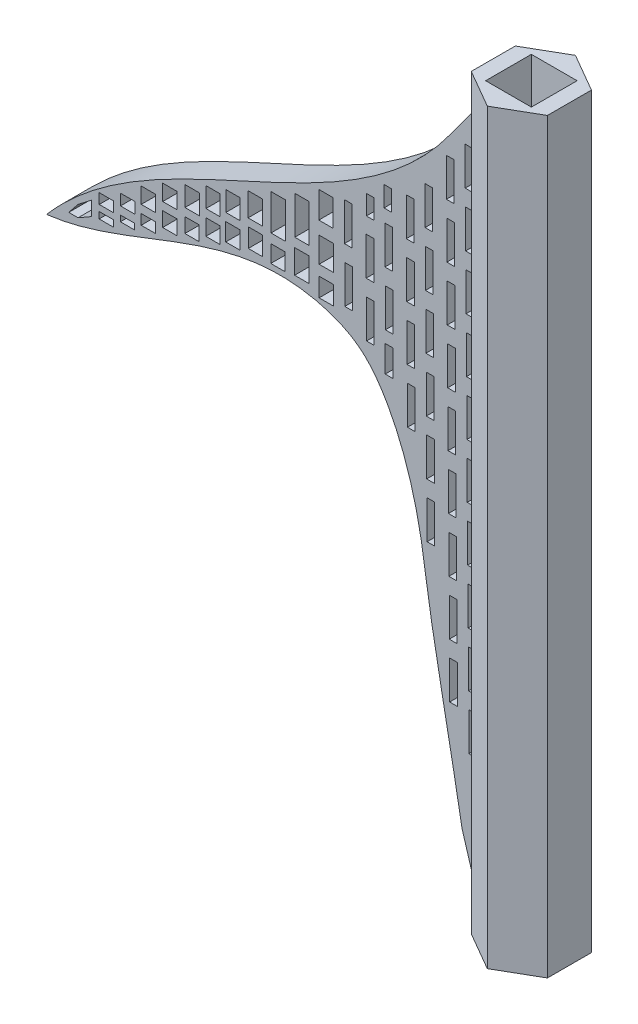
SolidWorks part; units mm, degrees
ref_plane "Front Plane" through (0, 0, 0) normal (0, 0, 1) x (1, 0, 0)
ref_plane "Top Plane" through (0, 0, 0) normal (0, 1, 0) x (1, 0, 0)
ref_plane "Right Plane" through (0, 0, 0) normal (1, 0, 0) x (0, 0, -1)
sketch "Sketch1" plane through (0, 0, 0) normal (0, 0, 1) x (1, 0, 0)
  line L0 (0.5851, 135.3104) -> (0.5851, 14.6604)
  line L1 (0.5851, 14.6604) -> (-3.4173, 27.924)
  line L2 (0.5851, 135.3104) -> (-5.3603, 127.1973)
  spline S0 degree 3 poles (-5.3603, 127.1973) (-22.25, 103.7542) (-54.2123, 103.4579) (-72.6613, 81.9767) knots 0 0 0 0 1 1 1 1
  spline S1 degree 3 poles (-72.6613, 81.9767) (-59.1241, 83.593) (-42.9036, 95.757) (-21.6318, 90.6459) (-14.6372, 82.9484) (-10.7236, 70.9466) (-8.6165, 54.5095) (-4.9898, 37.0221) (-3.4173, 27.924) knots 0 0 0 0 0.357139 0.42407 0.534017 0.754058 0.800656 1 1 1 1
  point P5 (-48.8145, 87.4527)
  point P8 (-54.1138, 87.6293)
  point P11 (-31.3269, 92.5753)
  point P13 (0, 0)
  point P15 (0, 0)
  point P17 (-5.3603, 24.0378)
  point P19 (-11.8961, 59.3664)
  point P20 (-3.4173, 27.924)
  point P21 (0, 0)
  point P22 (-9.5998, 62.1927)
  point P23 (-16.8421, 84.6264)
  point P24 (-23.9079, 90.8089)
extrude "Boss-Extrude1" add sketch "Sketch1" along normal blind 5.08 contours S0 S1 L1 L0 L2
sketch "Sketch2" plane through (0, 0, 5.08) normal (0, 0, 1) x (1, 0, 0)
  line L1 (-2.9091, 126.9995) -> (-1.6391, 126.9995)
  line L2 (-2.9091, 126.9995) -> (-2.9091, 120.6495)
  line L3 (-2.9091, 120.6495) -> (-1.6391, 120.6495)
  line L4 (-1.6391, 126.9995) -> (-1.6391, 120.6495)
  line L539 (-6.0375, 123.8245) -> (-6.0375, 117.4745)
  line L540 (-6.0375, 123.8245) -> (-4.7675, 123.8245)
  line L541 (-4.7675, 123.8245) -> (-4.7675, 117.4745)
  line L542 (-6.0375, 117.4745) -> (-4.7675, 117.4745)
  line L551 (-9.5949, 117.9664) -> (-8.3249, 117.9664)
  line L552 (-9.5949, 117.9664) -> (-9.5949, 111.6164)
  line L553 (-9.5949, 111.6164) -> (-8.3249, 111.6164)
  line L554 (-8.3249, 117.9664) -> (-8.3249, 111.6164)
  line L555 (-12.7232, 114.7914) -> (-12.7232, 108.4414)
  line L556 (-12.7232, 114.7914) -> (-11.4532, 114.7914)
  line L557 (-11.4532, 114.7914) -> (-11.4532, 108.4414)
  line L558 (-12.7232, 108.4414) -> (-11.4532, 108.4414)
  line L559 (-9.5272, 108.9333) -> (-8.2572, 108.9333)
  line L560 (-9.5272, 108.9333) -> (-9.5272, 102.5833)
  line L561 (-9.5272, 102.5833) -> (-8.2572, 102.5833)
  line L562 (-8.2572, 108.9333) -> (-8.2572, 102.5833)
  line L563 (-12.6556, 105.7583) -> (-12.6556, 99.4083)
  line L564 (-12.6556, 105.7583) -> (-11.3856, 105.7583)
  line L565 (-11.3856, 105.7583) -> (-11.3856, 99.4083)
  line L566 (-12.6556, 99.4083) -> (-11.3856, 99.4083)
  line L567 (-9.4596, 99.9002) -> (-8.1896, 99.9002)
  line L568 (-9.4596, 99.9002) -> (-9.4596, 93.5502)
  line L569 (-9.4596, 93.5502) -> (-8.1896, 93.5502)
  line L570 (-8.1896, 99.9002) -> (-8.1896, 93.5502)
  line L571 (-12.588, 96.7252) -> (-12.588, 90.3752)
  line L572 (-12.588, 96.7252) -> (-11.318, 96.7252)
  line L573 (-11.318, 96.7252) -> (-11.318, 90.3752)
  line L574 (-12.588, 90.3752) -> (-11.318, 90.3752)
  line L575 (-9.392, 90.8671) -> (-8.122, 90.8671)
  line L576 (-9.392, 90.8671) -> (-9.392, 84.5171)
  line L577 (-9.392, 84.5171) -> (-8.122, 84.5171)
  line L578 (-8.122, 90.8671) -> (-8.122, 84.5171)
  line L579 (-12.5203, 87.6921) -> (-12.5203, 81.3421)
  line L580 (-12.5203, 87.6921) -> (-11.2503, 87.6921)
  line L581 (-11.2503, 87.6921) -> (-11.2503, 81.3421)
  line L582 (-12.5203, 81.3421) -> (-11.2503, 81.3421)
  line L583 (-9.3243, 81.834) -> (-8.0543, 81.834)
  line L584 (-9.3243, 81.834) -> (-9.3243, 75.484)
  line L585 (-9.3243, 75.484) -> (-8.0543, 75.484)
  line L586 (-8.0543, 81.834) -> (-8.0543, 75.484)
  line L591 (-9.2567, 72.8009) -> (-7.9867, 72.8009)
  line L592 (-9.2567, 72.8009) -> (-9.2567, 66.4509)
  line L593 (-9.2567, 66.4509) -> (-7.9867, 66.4509)
  line L594 (-7.9867, 72.8009) -> (-7.9867, 66.4509)
  line L639 (-2.8415, 117.9664) -> (-1.5715, 117.9664)
  line L640 (-2.8415, 117.9664) -> (-2.8415, 111.6164)
  line L641 (-2.8415, 111.6164) -> (-1.5715, 111.6164)
  line L642 (-1.5715, 117.9664) -> (-1.5715, 111.6164)
  line L643 (-5.9699, 114.7914) -> (-5.9699, 108.4414)
  line L644 (-5.9699, 114.7914) -> (-4.6999, 114.7914)
  line L645 (-4.6999, 114.7914) -> (-4.6999, 108.4414)
  line L646 (-5.9699, 108.4414) -> (-4.6999, 108.4414)
  line L647 (-2.7739, 108.9333) -> (-1.5039, 108.9333)
  line L648 (-2.7739, 108.9333) -> (-2.7739, 102.5833)
  line L649 (-2.7739, 102.5833) -> (-1.5039, 102.5833)
  line L650 (-1.5039, 108.9333) -> (-1.5039, 102.5833)
  line L651 (-5.9022, 105.7583) -> (-5.9022, 99.4083)
  line L652 (-5.9022, 105.7583) -> (-4.6322, 105.7583)
  line L653 (-4.6322, 105.7583) -> (-4.6322, 99.4083)
  line L654 (-5.9022, 99.4083) -> (-4.6322, 99.4083)
  line L655 (-2.7062, 99.9002) -> (-1.4362, 99.9002)
  line L656 (-2.7062, 99.9002) -> (-2.7062, 93.5502)
  line L657 (-2.7062, 93.5502) -> (-1.4362, 93.5502)
  line L658 (-1.4362, 99.9002) -> (-1.4362, 93.5502)
  line L659 (-5.8346, 96.7252) -> (-5.8346, 90.3752)
  line L660 (-5.8346, 96.7252) -> (-4.5646, 96.7252)
  line L661 (-4.5646, 96.7252) -> (-4.5646, 90.3752)
  line L662 (-5.8346, 90.3752) -> (-4.5646, 90.3752)
  line L663 (-2.6386, 90.8671) -> (-1.3686, 90.8671)
  line L664 (-2.6386, 90.8671) -> (-2.6386, 84.5171)
  line L665 (-2.6386, 84.5171) -> (-1.3686, 84.5171)
  line L666 (-1.3686, 90.8671) -> (-1.3686, 84.5171)
  line L667 (-5.767, 87.6921) -> (-5.767, 81.3421)
  line L668 (-5.767, 87.6921) -> (-4.497, 87.6921)
  line L669 (-4.497, 87.6921) -> (-4.497, 81.3421)
  line L670 (-5.767, 81.3421) -> (-4.497, 81.3421)
  line L671 (-2.571, 81.834) -> (-1.301, 81.834)
  line L672 (-2.571, 81.834) -> (-2.571, 75.484)
  line L673 (-2.571, 75.484) -> (-1.301, 75.484)
  line L674 (-1.301, 81.834) -> (-1.301, 75.484)
  line L675 (-5.6993, 78.659) -> (-5.6993, 72.309)
  line L676 (-5.6993, 78.659) -> (-4.4293, 78.659)
  line L677 (-4.4293, 78.659) -> (-4.4293, 72.309)
  line L678 (-5.6993, 72.309) -> (-4.4293, 72.309)
  line L679 (-2.5033, 72.8009) -> (-1.2333, 72.8009)
  line L680 (-2.5033, 72.8009) -> (-2.5033, 66.4509)
  line L681 (-2.5033, 66.4509) -> (-1.2333, 66.4509)
  line L682 (-1.2333, 72.8009) -> (-1.2333, 66.4509)
  line L683 (-5.6317, 69.6259) -> (-5.6317, 63.2759)
  line L684 (-5.6317, 69.6259) -> (-4.3617, 69.6259)
  line L685 (-4.3617, 69.6259) -> (-4.3617, 63.2759)
  line L686 (-5.6317, 63.2759) -> (-4.3617, 63.2759)
  line L687 (-2.4357, 63.7678) -> (-1.1657, 63.7678)
  line L688 (-2.4357, 63.7678) -> (-2.4357, 57.4178)
  line L689 (-2.4357, 57.4178) -> (-1.1657, 57.4178)
  line L690 (-1.1657, 63.7678) -> (-1.1657, 57.4178)
  line L691 (-5.5641, 60.5928) -> (-5.5641, 54.2428)
  line L692 (-5.5641, 60.5928) -> (-4.2941, 60.5928)
  line L693 (-4.2941, 60.5928) -> (-4.2941, 54.2428)
  line L694 (-5.5641, 54.2428) -> (-4.2941, 54.2428)
  line L695 (-2.3681, 54.7347) -> (-1.0981, 54.7347)
  line L696 (-2.3681, 54.7347) -> (-2.3681, 48.3847)
  line L697 (-2.3681, 48.3847) -> (-1.0981, 48.3847)
  line L698 (-1.0981, 54.7347) -> (-1.0981, 48.3847)
  line L699 (-5.4964, 51.5597) -> (-5.4964, 45.2097)
  line L700 (-5.4964, 51.5597) -> (-4.2264, 51.5597)
  line L701 (-4.2264, 51.5597) -> (-4.2264, 45.2097)
  line L702 (-5.4964, 45.2097) -> (-4.2264, 45.2097)
  line L703 (-2.3005, 45.7016) -> (-1.0305, 45.7016)
  line L704 (-2.3005, 45.7016) -> (-2.3005, 39.3516)
  line L705 (-2.3005, 39.3516) -> (-1.0305, 39.3516)
  line L706 (-1.0305, 45.7016) -> (-1.0305, 39.3516)
  line L711 (-2.2328, 36.6685) -> (-0.9628, 36.6685)
  line L712 (-2.2328, 36.6685) -> (-2.2328, 30.3185)
  line L713 (-2.2328, 30.3185) -> (-0.9628, 30.3185)
  line L714 (-0.9628, 36.6685) -> (-0.9628, 30.3185)
  line L1047 (-16.2806, 108.9333) -> (-15.0106, 108.9333)
  line L1048 (-16.2806, 108.9333) -> (-16.2806, 102.5833)
  line L1049 (-16.2806, 102.5833) -> (-15.0106, 102.5833)
  line L1050 (-15.0106, 108.9333) -> (-15.0106, 102.5833)
  line L1051 (-19.4089, 105.7583) -> (-19.4089, 99.4083)
  line L1052 (-19.4089, 105.7583) -> (-18.1389, 105.7583)
  line L1053 (-18.1389, 105.7583) -> (-18.1389, 99.4083)
  line L1054 (-19.4089, 99.4083) -> (-18.1389, 99.4083)
  line L1055 (-23.0339, 108.9333) -> (-21.7639, 108.9333)
  line L1056 (-23.0339, 108.9333) -> (-23.0339, 102.5833)
  line L1057 (-23.0339, 102.5833) -> (-21.7639, 102.5833)
  line L1058 (-21.7639, 108.9333) -> (-21.7639, 102.5833)
  line L1111 (-16.213, 99.9002) -> (-14.943, 99.9002)
  line L1112 (-16.213, 99.9002) -> (-16.213, 93.5502)
  line L1113 (-16.213, 93.5502) -> (-14.943, 93.5502)
  line L1114 (-14.943, 99.9002) -> (-14.943, 93.5502)
  line L1115 (-19.3413, 96.7252) -> (-19.3413, 90.3752)
  line L1116 (-19.3413, 96.7252) -> (-18.0713, 96.7252)
  line L1117 (-18.0713, 96.7252) -> (-18.0713, 90.3752)
  line L1118 (-19.3413, 90.3752) -> (-18.0713, 90.3752)
  line L1119 (-22.9663, 99.9002) -> (-21.6963, 99.9002)
  line L1120 (-22.9663, 99.9002) -> (-22.9663, 93.5502)
  line L1121 (-22.9663, 93.5502) -> (-21.6963, 93.5502)
  line L1122 (-21.6963, 99.9002) -> (-21.6963, 93.5502)
  line L1687 (-12.1145, 33.4935) -> (-12.1145, 27.1435) [skipped]
  line L1688 (-12.0469, 24.4604) -> (-12.0469, 18.1104) [skipped]
  line L1689 (-16.0101, 66.4509) -> (-14.7401, 66.4509) [skipped]
  line L1690 (-19.1384, 63.2759) -> (-17.8684, 63.2759) [skipped]
  line L1691 (-22.7634, 66.4509) -> (-21.4934, 66.4509) [skipped]
  line L1692 (-25.8918, 63.2759) -> (-24.6218, 63.2759) [skipped]
  line L1693 (-29.5168, 66.4509) -> (-28.2468, 66.4509) [skipped]
  line L1694 (-32.6451, 63.2759) -> (-31.3751, 63.2759) [skipped]
  line L1695 (-36.2701, 66.4509) -> (-35.0001, 66.4509) [skipped]
  line L1696 (-39.3985, 63.2759) -> (-38.1285, 63.2759) [skipped]
  line L1697 (-43.0235, 66.4509) -> (-41.7535, 66.4509) [skipped]
  line L1698 (-46.1519, 63.2759) -> (-44.8819, 63.2759) [skipped]
  line L1699 (-49.7769, 66.4509) -> (-48.5069, 66.4509) [skipped]
  line L1700 (-52.9052, 63.2759) -> (-51.6352, 63.2759) [skipped]
  line L1701 (-56.5302, 66.4509) -> (-55.2602, 66.4509) [skipped]
  line L1702 (-59.6586, 63.2759) -> (-58.3886, 63.2759) [skipped]
  line L1703 (-63.2836, 66.4509) -> (-62.0136, 66.4509) [skipped]
  line L1704 (-66.4119, 63.2759) -> (-65.1419, 63.2759) [skipped]
  line L1705 (-15.9424, 63.7678) -> (-14.6724, 63.7678) [skipped]
  line L1706 (-15.9424, 63.7678) -> (-15.9424, 57.4178) [skipped]
  line L1707 (-15.9424, 57.4178) -> (-14.6724, 57.4178) [skipped]
  line L1708 (-14.6724, 63.7678) -> (-14.6724, 57.4178) [skipped]
  line L1709 (-19.0708, 60.5928) -> (-19.0708, 54.2428) [skipped]
  line L1710 (-19.0708, 60.5928) -> (-17.8008, 60.5928) [skipped]
  line L1711 (-17.8008, 60.5928) -> (-17.8008, 54.2428) [skipped]
  line L1712 (-19.0708, 54.2428) -> (-17.8008, 54.2428) [skipped]
  line L1713 (-22.6958, 63.7678) -> (-21.4258, 63.7678) [skipped]
  line L1714 (-22.6958, 63.7678) -> (-22.6958, 57.4178) [skipped]
  line L1715 (-22.6958, 57.4178) -> (-21.4258, 57.4178) [skipped]
  line L1716 (-21.4258, 63.7678) -> (-21.4258, 57.4178) [skipped]
  line L1717 (-25.8241, 60.5928) -> (-25.8241, 54.2428) [skipped]
  line L1718 (-25.8241, 60.5928) -> (-24.5541, 60.5928) [skipped]
  line L1719 (-24.5541, 60.5928) -> (-24.5541, 54.2428) [skipped]
  line L1720 (-25.8241, 54.2428) -> (-24.5541, 54.2428) [skipped]
  line L1721 (-29.4491, 63.7678) -> (-28.1791, 63.7678) [skipped]
  line L1722 (-29.4491, 63.7678) -> (-29.4491, 57.4178) [skipped]
  line L1723 (-29.4491, 57.4178) -> (-28.1791, 57.4178) [skipped]
  line L1724 (-28.1791, 63.7678) -> (-28.1791, 57.4178) [skipped]
  line L1725 (-32.5775, 60.5928) -> (-32.5775, 54.2428) [skipped]
  line L1726 (-32.5775, 60.5928) -> (-31.3075, 60.5928) [skipped]
  line L1727 (-31.3075, 60.5928) -> (-31.3075, 54.2428) [skipped]
  line L1728 (-32.5775, 54.2428) -> (-31.3075, 54.2428) [skipped]
  line L1729 (-36.2025, 63.7678) -> (-34.9325, 63.7678) [skipped]
  line L1730 (-36.2025, 63.7678) -> (-36.2025, 57.4178) [skipped]
  line L1731 (-36.2025, 57.4178) -> (-34.9325, 57.4178) [skipped]
  line L1732 (-34.9325, 63.7678) -> (-34.9325, 57.4178) [skipped]
  line L1733 (-39.3309, 60.5928) -> (-39.3309, 54.2428) [skipped]
  line L1734 (-39.3309, 60.5928) -> (-38.0609, 60.5928) [skipped]
  line L1735 (-38.0609, 60.5928) -> (-38.0609, 54.2428) [skipped]
  line L1736 (-39.3309, 54.2428) -> (-38.0609, 54.2428) [skipped]
  line L1737 (-42.9559, 63.7678) -> (-41.6859, 63.7678) [skipped]
  line L1738 (-42.9559, 63.7678) -> (-42.9559, 57.4178) [skipped]
  line L1739 (-42.9559, 57.4178) -> (-41.6859, 57.4178) [skipped]
  line L1740 (-41.6859, 63.7678) -> (-41.6859, 57.4178) [skipped]
  line L1741 (-46.0842, 60.5928) -> (-46.0842, 54.2428) [skipped]
  line L1742 (-46.0842, 60.5928) -> (-44.8142, 60.5928) [skipped]
  line L1743 (-44.8142, 60.5928) -> (-44.8142, 54.2428) [skipped]
  line L1744 (-46.0842, 54.2428) -> (-44.8142, 54.2428) [skipped]
  line L1745 (-49.7092, 63.7678) -> (-48.4392, 63.7678) [skipped]
  line L1746 (-49.7092, 63.7678) -> (-49.7092, 57.4178) [skipped]
  line L1747 (-49.7092, 57.4178) -> (-48.4392, 57.4178) [skipped]
  line L1748 (-48.4392, 63.7678) -> (-48.4392, 57.4178) [skipped]
  line L1749 (-52.8376, 60.5928) -> (-52.8376, 54.2428) [skipped]
  line L1750 (-52.8376, 60.5928) -> (-51.5676, 60.5928) [skipped]
  line L1751 (-51.5676, 60.5928) -> (-51.5676, 54.2428) [skipped]
  line L1752 (-52.8376, 54.2428) -> (-51.5676, 54.2428) [skipped]
  line L1753 (-56.4626, 63.7678) -> (-55.1926, 63.7678) [skipped]
  line L1754 (-56.4626, 63.7678) -> (-56.4626, 57.4178) [skipped]
  line L1755 (-56.4626, 57.4178) -> (-55.1926, 57.4178) [skipped]
  line L1756 (-55.1926, 63.7678) -> (-55.1926, 57.4178) [skipped]
  line L1757 (-59.5909, 60.5928) -> (-59.5909, 54.2428) [skipped]
  line L1758 (-59.5909, 60.5928) -> (-58.3209, 60.5928) [skipped]
  line L1759 (-58.3209, 60.5928) -> (-58.3209, 54.2428) [skipped]
  line L1760 (-59.5909, 54.2428) -> (-58.3209, 54.2428) [skipped]
  line L1761 (-63.2159, 63.7678) -> (-61.9459, 63.7678) [skipped]
  line L1762 (-63.2159, 63.7678) -> (-63.2159, 57.4178) [skipped]
  line L1763 (-63.2159, 57.4178) -> (-61.9459, 57.4178) [skipped]
  line L1764 (-61.9459, 63.7678) -> (-61.9459, 57.4178) [skipped]
  line L1765 (-66.3443, 60.5928) -> (-66.3443, 54.2428) [skipped]
  line L1766 (-66.3443, 60.5928) -> (-65.0743, 60.5928) [skipped]
  line L1767 (-65.0743, 60.5928) -> (-65.0743, 54.2428) [skipped]
  line L1768 (-66.3443, 54.2428) -> (-65.0743, 54.2428) [skipped]
  line L1769 (-15.8748, 54.7347) -> (-14.6048, 54.7347) [skipped]
  line L1770 (-15.8748, 54.7347) -> (-15.8748, 48.3847) [skipped]
  line L1771 (-15.8748, 48.3847) -> (-14.6048, 48.3847) [skipped]
  line L1772 (-14.6048, 54.7347) -> (-14.6048, 48.3847) [skipped]
  line L1773 (-19.0032, 51.5597) -> (-19.0032, 45.2097) [skipped]
  line L1774 (-19.0032, 51.5597) -> (-17.7332, 51.5597) [skipped]
  line L1775 (-17.7332, 51.5597) -> (-17.7332, 45.2097) [skipped]
  line L1776 (-19.0032, 45.2097) -> (-17.7332, 45.2097) [skipped]
  line L1777 (-22.6282, 54.7347) -> (-21.3582, 54.7347) [skipped]
  line L1778 (-22.6282, 54.7347) -> (-22.6282, 48.3847) [skipped]
  line L1779 (-22.6282, 48.3847) -> (-21.3582, 48.3847) [skipped]
  line L1780 (-21.3582, 54.7347) -> (-21.3582, 48.3847) [skipped]
  line L1781 (-25.7565, 51.5597) -> (-25.7565, 45.2097) [skipped]
  line L1782 (-25.7565, 51.5597) -> (-24.4865, 51.5597) [skipped]
  line L1783 (-24.4865, 51.5597) -> (-24.4865, 45.2097) [skipped]
  line L1784 (-25.7565, 45.2097) -> (-24.4865, 45.2097) [skipped]
  line L1785 (-29.3815, 54.7347) -> (-28.1115, 54.7347) [skipped]
  line L1786 (-29.3815, 54.7347) -> (-29.3815, 48.3847) [skipped]
  line L1787 (-29.3815, 48.3847) -> (-28.1115, 48.3847) [skipped]
  line L1788 (-28.1115, 54.7347) -> (-28.1115, 48.3847) [skipped]
  line L1789 (-32.5099, 51.5597) -> (-32.5099, 45.2097) [skipped]
  line L1790 (-32.5099, 51.5597) -> (-31.2399, 51.5597) [skipped]
  line L1791 (-31.2399, 51.5597) -> (-31.2399, 45.2097) [skipped]
  line L1792 (-32.5099, 45.2097) -> (-31.2399, 45.2097) [skipped]
  line L1793 (-36.1349, 54.7347) -> (-34.8649, 54.7347) [skipped]
  line L1794 (-36.1349, 54.7347) -> (-36.1349, 48.3847) [skipped]
  line L1795 (-36.1349, 48.3847) -> (-34.8649, 48.3847) [skipped]
  line L1796 (-34.8649, 54.7347) -> (-34.8649, 48.3847) [skipped]
  line L1797 (-39.2632, 51.5597) -> (-39.2632, 45.2097) [skipped]
  line L1798 (-39.2632, 51.5597) -> (-37.9932, 51.5597) [skipped]
  line L1799 (-37.9932, 51.5597) -> (-37.9932, 45.2097) [skipped]
  line L1800 (-39.2632, 45.2097) -> (-37.9932, 45.2097) [skipped]
  line L1801 (-42.8882, 54.7347) -> (-41.6182, 54.7347) [skipped]
  line L1802 (-42.8882, 54.7347) -> (-42.8882, 48.3847) [skipped]
  line L1803 (-42.8882, 48.3847) -> (-41.6182, 48.3847) [skipped]
  line L1804 (-41.6182, 54.7347) -> (-41.6182, 48.3847) [skipped]
  line L1805 (-46.0166, 51.5597) -> (-46.0166, 45.2097) [skipped]
  line L1806 (-46.0166, 51.5597) -> (-44.7466, 51.5597) [skipped]
  line L1807 (-44.7466, 51.5597) -> (-44.7466, 45.2097) [skipped]
  line L1808 (-46.0166, 45.2097) -> (-44.7466, 45.2097) [skipped]
  line L1809 (-49.6416, 54.7347) -> (-48.3716, 54.7347) [skipped]
  line L1810 (-49.6416, 54.7347) -> (-49.6416, 48.3847) [skipped]
  line L1811 (-49.6416, 48.3847) -> (-48.3716, 48.3847) [skipped]
  line L1812 (-48.3716, 54.7347) -> (-48.3716, 48.3847) [skipped]
  line L1813 (-52.7699, 51.5597) -> (-52.7699, 45.2097) [skipped]
  line L1814 (-52.7699, 51.5597) -> (-51.4999, 51.5597) [skipped]
  line L1815 (-51.4999, 51.5597) -> (-51.4999, 45.2097) [skipped]
  line L1816 (-52.7699, 45.2097) -> (-51.4999, 45.2097) [skipped]
  line L1817 (-56.395, 54.7347) -> (-55.125, 54.7347) [skipped]
  line L1818 (-56.395, 54.7347) -> (-56.395, 48.3847) [skipped]
  line L1819 (-56.395, 48.3847) -> (-55.125, 48.3847) [skipped]
  line L1820 (-55.125, 54.7347) -> (-55.125, 48.3847) [skipped]
  line L1821 (-59.5233, 51.5597) -> (-59.5233, 45.2097) [skipped]
  line L1822 (-59.5233, 51.5597) -> (-58.2533, 51.5597) [skipped]
  line L1823 (-58.2533, 51.5597) -> (-58.2533, 45.2097) [skipped]
  line L1824 (-59.5233, 45.2097) -> (-58.2533, 45.2097) [skipped]
  line L1825 (-63.1483, 54.7347) -> (-61.8783, 54.7347) [skipped]
  line L1826 (-63.1483, 54.7347) -> (-63.1483, 48.3847) [skipped]
  line L1827 (-63.1483, 48.3847) -> (-61.8783, 48.3847) [skipped]
  line L1828 (-61.8783, 54.7347) -> (-61.8783, 48.3847) [skipped]
  line L1829 (-66.2767, 51.5597) -> (-66.2767, 45.2097) [skipped]
  line L1830 (-66.2767, 51.5597) -> (-65.0067, 51.5597) [skipped]
  line L1831 (-65.0067, 51.5597) -> (-65.0067, 45.2097) [skipped]
  line L1832 (-66.2767, 45.2097) -> (-65.0067, 45.2097) [skipped]
  line L1833 (-15.8072, 45.7016) -> (-14.5372, 45.7016) [skipped]
  line L1834 (-15.8072, 45.7016) -> (-15.8072, 39.3516) [skipped]
  line L1835 (-15.8072, 39.3516) -> (-14.5372, 39.3516) [skipped]
  line L1836 (-14.5372, 45.7016) -> (-14.5372, 39.3516) [skipped]
  line L1837 (-18.9355, 42.5266) -> (-18.9355, 36.1766) [skipped]
  line L1838 (-18.9355, 42.5266) -> (-17.6655, 42.5266) [skipped]
  line L1839 (-17.6655, 42.5266) -> (-17.6655, 36.1766) [skipped]
  line L1840 (-18.9355, 36.1766) -> (-17.6655, 36.1766) [skipped]
  line L1841 (-22.5605, 45.7016) -> (-21.2905, 45.7016) [skipped]
  line L1842 (-22.5605, 45.7016) -> (-22.5605, 39.3516) [skipped]
  line L1843 (-22.5605, 39.3516) -> (-21.2905, 39.3516) [skipped]
  line L1844 (-21.2905, 45.7016) -> (-21.2905, 39.3516) [skipped]
  line L1845 (-25.6889, 42.5266) -> (-25.6889, 36.1766) [skipped]
  line L1846 (-25.6889, 42.5266) -> (-24.4189, 42.5266) [skipped]
  line L1847 (-24.4189, 42.5266) -> (-24.4189, 36.1766) [skipped]
  line L1848 (-25.6889, 36.1766) -> (-24.4189, 36.1766) [skipped]
  line L1849 (-29.3139, 45.7016) -> (-28.0439, 45.7016) [skipped]
  line L1850 (-29.3139, 45.7016) -> (-29.3139, 39.3516) [skipped]
  line L1851 (-29.3139, 39.3516) -> (-28.0439, 39.3516) [skipped]
  line L1852 (-28.0439, 45.7016) -> (-28.0439, 39.3516) [skipped]
  line L1853 (-32.4422, 42.5266) -> (-32.4422, 36.1766) [skipped]
  line L1854 (-32.4422, 42.5266) -> (-31.1722, 42.5266) [skipped]
  line L1855 (-31.1722, 42.5266) -> (-31.1722, 36.1766) [skipped]
  line L1856 (-32.4422, 36.1766) -> (-31.1722, 36.1766) [skipped]
  line L1857 (-36.0672, 45.7016) -> (-34.7972, 45.7016) [skipped]
  line L1858 (-36.0672, 45.7016) -> (-36.0672, 39.3516) [skipped]
  line L1859 (-36.0672, 39.3516) -> (-34.7972, 39.3516) [skipped]
  line L1860 (-34.7972, 45.7016) -> (-34.7972, 39.3516) [skipped]
  line L1861 (-39.1956, 42.5266) -> (-39.1956, 36.1766) [skipped]
  line L1862 (-39.1956, 42.5266) -> (-37.9256, 42.5266) [skipped]
  line L1863 (-37.9256, 42.5266) -> (-37.9256, 36.1766) [skipped]
  line L1864 (-39.1956, 36.1766) -> (-37.9256, 36.1766) [skipped]
  line L1865 (-42.8206, 45.7016) -> (-41.5506, 45.7016) [skipped]
  line L1866 (-42.8206, 45.7016) -> (-42.8206, 39.3516) [skipped]
  line L1867 (-42.8206, 39.3516) -> (-41.5506, 39.3516) [skipped]
  line L1868 (-41.5506, 45.7016) -> (-41.5506, 39.3516) [skipped]
  line L1869 (-45.949, 42.5266) -> (-45.949, 36.1766) [skipped]
  line L1870 (-45.949, 42.5266) -> (-44.679, 42.5266) [skipped]
  line L1871 (-44.679, 42.5266) -> (-44.679, 36.1766) [skipped]
  line L1872 (-45.949, 36.1766) -> (-44.679, 36.1766) [skipped]
  line L1873 (-49.574, 45.7016) -> (-48.304, 45.7016) [skipped]
  line L1874 (-49.574, 45.7016) -> (-49.574, 39.3516) [skipped]
  line L1875 (-49.574, 39.3516) -> (-48.304, 39.3516) [skipped]
  line L1876 (-48.304, 45.7016) -> (-48.304, 39.3516) [skipped]
  line L1877 (-52.7023, 42.5266) -> (-52.7023, 36.1766) [skipped]
  line L1878 (-52.7023, 42.5266) -> (-51.4323, 42.5266) [skipped]
  line L1879 (-51.4323, 42.5266) -> (-51.4323, 36.1766) [skipped]
  line L1880 (-52.7023, 36.1766) -> (-51.4323, 36.1766) [skipped]
  line L1881 (-56.3273, 45.7016) -> (-55.0573, 45.7016) [skipped]
  line L1882 (-56.3273, 45.7016) -> (-56.3273, 39.3516) [skipped]
  line L1883 (-56.3273, 39.3516) -> (-55.0573, 39.3516) [skipped]
  line L1884 (-55.0573, 45.7016) -> (-55.0573, 39.3516) [skipped]
  line L1885 (-59.4557, 42.5266) -> (-59.4557, 36.1766) [skipped]
  line L1886 (-59.4557, 42.5266) -> (-58.1857, 42.5266) [skipped]
  line L1887 (-58.1857, 42.5266) -> (-58.1857, 36.1766) [skipped]
  line L1888 (-59.4557, 36.1766) -> (-58.1857, 36.1766) [skipped]
  line L1889 (-63.0807, 45.7016) -> (-61.8107, 45.7016) [skipped]
  line L1890 (-63.0807, 45.7016) -> (-63.0807, 39.3516) [skipped]
  line L1891 (-63.0807, 39.3516) -> (-61.8107, 39.3516) [skipped]
  line L1892 (-61.8107, 45.7016) -> (-61.8107, 39.3516) [skipped]
  line L1893 (-66.209, 42.5266) -> (-66.209, 36.1766) [skipped]
  line L1894 (-66.209, 42.5266) -> (-64.939, 42.5266) [skipped]
  line L1895 (-64.939, 42.5266) -> (-64.939, 36.1766) [skipped]
  line L1896 (-66.209, 36.1766) -> (-64.939, 36.1766) [skipped]
  line L1897 (-15.7395, 36.6685) -> (-14.4695, 36.6685) [skipped]
  line L1898 (-15.7395, 36.6685) -> (-15.7395, 30.3185) [skipped]
  line L1899 (-15.7395, 30.3185) -> (-14.4695, 30.3185) [skipped]
  line L1900 (-14.4695, 36.6685) -> (-14.4695, 30.3185) [skipped]
  line L1901 (-18.8679, 33.4935) -> (-18.8679, 27.1435) [skipped]
  line L1902 (-18.8679, 33.4935) -> (-17.5979, 33.4935) [skipped]
  line L1903 (-17.5979, 33.4935) -> (-17.5979, 27.1435) [skipped]
  line L1904 (-18.8679, 27.1435) -> (-17.5979, 27.1435) [skipped]
  line L1905 (-22.4929, 36.6685) -> (-21.2229, 36.6685) [skipped]
  line L1906 (-22.4929, 36.6685) -> (-22.4929, 30.3185) [skipped]
  line L1907 (-22.4929, 30.3185) -> (-21.2229, 30.3185) [skipped]
  line L1908 (-21.2229, 36.6685) -> (-21.2229, 30.3185) [skipped]
  line L1909 (-25.6213, 33.4935) -> (-25.6213, 27.1435) [skipped]
  line L1910 (-25.6213, 33.4935) -> (-24.3513, 33.4935) [skipped]
  line L1911 (-24.3513, 33.4935) -> (-24.3513, 27.1435) [skipped]
  line L1912 (-25.6213, 27.1435) -> (-24.3513, 27.1435) [skipped]
  line L1913 (-29.2463, 36.6685) -> (-27.9763, 36.6685) [skipped]
  line L1914 (-29.2463, 36.6685) -> (-29.2463, 30.3185) [skipped]
  line L1915 (-29.2463, 30.3185) -> (-27.9763, 30.3185) [skipped]
  line L1916 (-27.9763, 36.6685) -> (-27.9763, 30.3185) [skipped]
  line L1917 (-32.3746, 33.4935) -> (-32.3746, 27.1435) [skipped]
  line L1918 (-32.3746, 33.4935) -> (-31.1046, 33.4935) [skipped]
  line L1919 (-31.1046, 33.4935) -> (-31.1046, 27.1435) [skipped]
  line L1920 (-32.3746, 27.1435) -> (-31.1046, 27.1435) [skipped]
  line L1921 (-35.9996, 36.6685) -> (-34.7296, 36.6685) [skipped]
  line L1922 (-35.9996, 36.6685) -> (-35.9996, 30.3185) [skipped]
  line L1923 (-35.9996, 30.3185) -> (-34.7296, 30.3185) [skipped]
  line L1924 (-34.7296, 36.6685) -> (-34.7296, 30.3185) [skipped]
  line L1925 (-39.128, 33.4935) -> (-39.128, 27.1435) [skipped]
  line L1926 (-39.128, 33.4935) -> (-37.858, 33.4935) [skipped]
  line L1927 (-37.858, 33.4935) -> (-37.858, 27.1435) [skipped]
  line L1928 (-39.128, 27.1435) -> (-37.858, 27.1435) [skipped]
  line L1929 (-42.753, 36.6685) -> (-41.483, 36.6685) [skipped]
  line L1930 (-42.753, 36.6685) -> (-42.753, 30.3185) [skipped]
  line L1931 (-42.753, 30.3185) -> (-41.483, 30.3185) [skipped]
  line L1932 (-41.483, 36.6685) -> (-41.483, 30.3185) [skipped]
  line L1933 (-45.8813, 33.4935) -> (-45.8813, 27.1435) [skipped]
  line L1934 (-45.8813, 33.4935) -> (-44.6113, 33.4935) [skipped]
  line L1935 (-44.6113, 33.4935) -> (-44.6113, 27.1435) [skipped]
  line L1936 (-45.8813, 27.1435) -> (-44.6113, 27.1435) [skipped]
  line L1937 (-49.5063, 36.6685) -> (-48.2363, 36.6685) [skipped]
  line L1938 (-49.5063, 36.6685) -> (-49.5063, 30.3185) [skipped]
  line L1939 (-49.5063, 30.3185) -> (-48.2363, 30.3185) [skipped]
  line L1940 (-48.2363, 36.6685) -> (-48.2363, 30.3185) [skipped]
  line L1941 (-52.6347, 33.4935) -> (-52.6347, 27.1435) [skipped]
  line L1942 (-52.6347, 33.4935) -> (-51.3647, 33.4935) [skipped]
  line L1943 (-51.3647, 33.4935) -> (-51.3647, 27.1435) [skipped]
  line L1944 (-52.6347, 27.1435) -> (-51.3647, 27.1435) [skipped]
  line L1945 (-56.2597, 36.6685) -> (-54.9897, 36.6685) [skipped]
  line L1946 (-56.2597, 36.6685) -> (-56.2597, 30.3185) [skipped]
  line L1947 (-56.2597, 30.3185) -> (-54.9897, 30.3185) [skipped]
  line L1948 (-54.9897, 36.6685) -> (-54.9897, 30.3185) [skipped]
  line L1949 (-59.388, 33.4935) -> (-59.388, 27.1435) [skipped]
  line L1950 (-59.388, 33.4935) -> (-58.118, 33.4935) [skipped]
  line L1951 (-58.118, 33.4935) -> (-58.118, 27.1435) [skipped]
  line L1952 (-59.388, 27.1435) -> (-58.118, 27.1435) [skipped]
  line L1953 (-63.013, 36.6685) -> (-61.743, 36.6685) [skipped]
  line L1954 (-63.013, 36.6685) -> (-63.013, 30.3185) [skipped]
  line L1955 (-63.013, 30.3185) -> (-61.743, 30.3185) [skipped]
  line L1956 (-61.743, 36.6685) -> (-61.743, 30.3185) [skipped]
  line L1957 (-66.1414, 33.4935) -> (-66.1414, 27.1435) [skipped]
  line L1958 (-66.1414, 33.4935) -> (-64.8714, 33.4935) [skipped]
  line L1959 (-64.8714, 33.4935) -> (-64.8714, 27.1435) [skipped]
  line L1960 (-66.1414, 27.1435) -> (-64.8714, 27.1435) [skipped]
  line L1961 (-15.6719, 27.6354) -> (-14.4019, 27.6354) [skipped]
  line L1962 (-15.6719, 27.6354) -> (-15.6719, 21.2854) [skipped]
  line L1963 (-15.6719, 21.2854) -> (-14.4019, 21.2854) [skipped]
  line L1964 (-14.4019, 27.6354) -> (-14.4019, 21.2854) [skipped]
  line L1965 (-18.8003, 24.4604) -> (-18.8003, 18.1104) [skipped]
  line L1966 (-18.8003, 24.4604) -> (-17.5303, 24.4604) [skipped]
  line L1967 (-17.5303, 24.4604) -> (-17.5303, 18.1104) [skipped]
  line L1968 (-18.8003, 18.1104) -> (-17.5303, 18.1104) [skipped]
  line L1969 (-22.4253, 27.6354) -> (-21.1553, 27.6354) [skipped]
  line L1970 (-22.4253, 27.6354) -> (-22.4253, 21.2854) [skipped]
  line L1971 (-22.4253, 21.2854) -> (-21.1553, 21.2854) [skipped]
  line L1972 (-21.1553, 27.6354) -> (-21.1553, 21.2854) [skipped]
  line L1973 (-25.5536, 24.4604) -> (-25.5536, 18.1104) [skipped]
  line L1974 (-25.5536, 24.4604) -> (-24.2836, 24.4604) [skipped]
  line L1975 (-24.2836, 24.4604) -> (-24.2836, 18.1104) [skipped]
  line L1976 (-25.5536, 18.1104) -> (-24.2836, 18.1104) [skipped]
  line L1977 (-29.1786, 27.6354) -> (-27.9086, 27.6354) [skipped]
  line L1978 (-29.1786, 27.6354) -> (-29.1786, 21.2854) [skipped]
  line L1979 (-29.1786, 21.2854) -> (-27.9086, 21.2854) [skipped]
  line L1980 (-27.9086, 27.6354) -> (-27.9086, 21.2854) [skipped]
  line L1981 (-32.307, 24.4604) -> (-32.307, 18.1104) [skipped]
  line L1982 (-32.307, 24.4604) -> (-31.037, 24.4604) [skipped]
  line L1983 (-31.037, 24.4604) -> (-31.037, 18.1104) [skipped]
  line L1984 (-32.307, 18.1104) -> (-31.037, 18.1104) [skipped]
  line L1985 (-35.932, 27.6354) -> (-34.662, 27.6354) [skipped]
  line L1986 (-35.932, 27.6354) -> (-35.932, 21.2854) [skipped]
  line L1987 (-35.932, 21.2854) -> (-34.662, 21.2854) [skipped]
  line L1988 (-34.662, 27.6354) -> (-34.662, 21.2854) [skipped]
  line L1989 (-39.0603, 24.4604) -> (-39.0603, 18.1104) [skipped]
  line L1990 (-39.0603, 24.4604) -> (-37.7903, 24.4604) [skipped]
  line L1991 (-37.7903, 24.4604) -> (-37.7903, 18.1104) [skipped]
  line L1992 (-39.0603, 18.1104) -> (-37.7903, 18.1104) [skipped]
  line L1993 (-42.6853, 27.6354) -> (-41.4153, 27.6354) [skipped]
  line L1994 (-42.6853, 27.6354) -> (-42.6853, 21.2854) [skipped]
  line L1995 (-42.6853, 21.2854) -> (-41.4153, 21.2854) [skipped]
  line L1996 (-41.4153, 27.6354) -> (-41.4153, 21.2854) [skipped]
  line L1997 (-45.8137, 24.4604) -> (-45.8137, 18.1104) [skipped]
  line L1998 (-45.8137, 24.4604) -> (-44.5437, 24.4604) [skipped]
  line L1999 (-44.5437, 24.4604) -> (-44.5437, 18.1104) [skipped]
  line L2000 (-45.8137, 18.1104) -> (-44.5437, 18.1104) [skipped]
  line L2001 (-49.4387, 27.6354) -> (-48.1687, 27.6354) [skipped]
  line L2002 (-49.4387, 27.6354) -> (-49.4387, 21.2854) [skipped]
  line L2003 (-49.4387, 21.2854) -> (-48.1687, 21.2854) [skipped]
  line L2004 (-48.1687, 27.6354) -> (-48.1687, 21.2854) [skipped]
  line L2005 (-52.5671, 24.4604) -> (-52.5671, 18.1104) [skipped]
  line L2006 (-52.5671, 24.4604) -> (-51.2971, 24.4604) [skipped]
  line L2007 (-51.2971, 24.4604) -> (-51.2971, 18.1104) [skipped]
  line L2008 (-52.5671, 18.1104) -> (-51.2971, 18.1104) [skipped]
  line L2009 (-56.1921, 27.6354) -> (-54.9221, 27.6354) [skipped]
  line L2010 (-56.1921, 27.6354) -> (-56.1921, 21.2854) [skipped]
  line L2011 (-56.1921, 21.2854) -> (-54.9221, 21.2854) [skipped]
  line L2012 (-54.9221, 27.6354) -> (-54.9221, 21.2854) [skipped]
  line L2013 (-59.3204, 24.4604) -> (-59.3204, 18.1104) [skipped]
  line L2014 (-59.3204, 24.4604) -> (-58.0504, 24.4604) [skipped]
  line L2015 (-58.0504, 24.4604) -> (-58.0504, 18.1104) [skipped]
  line L2016 (-59.3204, 18.1104) -> (-58.0504, 18.1104) [skipped]
  line L2017 (-62.9454, 27.6354) -> (-61.6754, 27.6354) [skipped]
  line L2018 (-62.9454, 27.6354) -> (-62.9454, 21.2854) [skipped]
  line L2019 (-62.9454, 21.2854) -> (-61.6754, 21.2854) [skipped]
  line L2020 (-61.6754, 27.6354) -> (-61.6754, 21.2854) [skipped]
  line L2021 (-66.0738, 24.4604) -> (-66.0738, 18.1104) [skipped]
  line L2022 (-66.0738, 24.4604) -> (-64.8038, 24.4604) [skipped]
  line L2023 (-64.8038, 24.4604) -> (-64.8038, 18.1104) [skipped]
  line L2024 (-66.0738, 18.1104) -> (-64.8038, 18.1104) [skipped]
  line L2025 (-33.0509, 123.8245) -> (-33.0509, 117.4745) [skipped]
  line L2026 (-36.6759, 126.9995) -> (-35.4059, 126.9995) [skipped]
  line L2027 (-36.6759, 126.9995) -> (-36.6759, 120.6495) [skipped]
  line L2028 (-36.6759, 120.6495) -> (-35.4059, 120.6495) [skipped]
  line L2029 (-35.4059, 126.9995) -> (-35.4059, 120.6495) [skipped]
  line L2030 (-39.8043, 123.8245) -> (-39.8043, 117.4745) [skipped]
  line L2031 (-39.8043, 123.8245) -> (-38.5343, 123.8245) [skipped]
  line L2032 (-38.5343, 123.8245) -> (-38.5343, 117.4745) [skipped]
  line L2033 (-39.8043, 117.4745) -> (-38.5343, 117.4745) [skipped]
  line L2034 (-43.4293, 126.9995) -> (-42.1593, 126.9995) [skipped]
  line L2035 (-43.4293, 126.9995) -> (-43.4293, 120.6495) [skipped]
  line L2036 (-43.4293, 120.6495) -> (-42.1593, 120.6495) [skipped]
  line L2037 (-42.1593, 126.9995) -> (-42.1593, 120.6495) [skipped]
  line L2038 (-46.5576, 123.8245) -> (-46.5576, 117.4745) [skipped]
  line L2039 (-46.5576, 123.8245) -> (-45.2876, 123.8245) [skipped]
  line L2040 (-45.2876, 123.8245) -> (-45.2876, 117.4745) [skipped]
  line L2041 (-46.5576, 117.4745) -> (-45.2876, 117.4745) [skipped]
  line L2042 (-50.1826, 126.9995) -> (-48.9126, 126.9995) [skipped]
  line L2043 (-50.1826, 126.9995) -> (-50.1826, 120.6495) [skipped]
  line L2044 (-50.1826, 120.6495) -> (-48.9126, 120.6495) [skipped]
  line L2045 (-48.9126, 126.9995) -> (-48.9126, 120.6495) [skipped]
  line L2046 (-53.311, 123.8245) -> (-53.311, 117.4745) [skipped]
  line L2047 (-53.311, 123.8245) -> (-52.041, 123.8245) [skipped]
  line L2048 (-52.041, 123.8245) -> (-52.041, 117.4745) [skipped]
  line L2049 (-53.311, 117.4745) -> (-52.041, 117.4745) [skipped]
  line L2050 (-56.936, 126.9995) -> (-55.666, 126.9995) [skipped]
  line L2051 (-56.936, 126.9995) -> (-56.936, 120.6495) [skipped]
  line L2052 (-56.936, 120.6495) -> (-55.666, 120.6495) [skipped]
  line L2053 (-55.666, 126.9995) -> (-55.666, 120.6495) [skipped]
  line L2054 (-60.0644, 123.8245) -> (-60.0644, 117.4745) [skipped]
  line L2055 (-60.0644, 123.8245) -> (-58.7944, 123.8245) [skipped]
  line L2056 (-58.7944, 123.8245) -> (-58.7944, 117.4745) [skipped]
  line L2057 (-60.0644, 117.4745) -> (-58.7944, 117.4745) [skipped]
  line L2058 (-63.6894, 126.9995) -> (-62.4194, 126.9995) [skipped]
  line L2059 (-63.6894, 126.9995) -> (-63.6894, 120.6495) [skipped]
  line L2060 (-63.6894, 120.6495) -> (-62.4194, 120.6495) [skipped]
  line L2061 (-62.4194, 126.9995) -> (-62.4194, 120.6495) [skipped]
  line L2062 (-66.8177, 123.8245) -> (-66.8177, 117.4745) [skipped]
  line L2063 (-66.8177, 123.8245) -> (-65.5477, 123.8245) [skipped]
  line L2064 (-65.5477, 123.8245) -> (-65.5477, 117.4745) [skipped]
  line L2065 (-66.8177, 117.4745) -> (-65.5477, 117.4745) [skipped]
  line L2066 (-36.6083, 117.9664) -> (-35.3383, 117.9664) [skipped]
  line L2067 (-36.6083, 117.9664) -> (-36.6083, 111.6164) [skipped]
  line L2068 (-36.6083, 111.6164) -> (-35.3383, 111.6164) [skipped]
  line L2069 (-35.3383, 117.9664) -> (-35.3383, 111.6164) [skipped]
  line L2070 (-39.7367, 114.7914) -> (-38.4667, 114.7914) [skipped]
  line L2071 (-43.3617, 117.9664) -> (-42.0917, 117.9664) [skipped]
  line L2072 (-43.3617, 117.9664) -> (-43.3617, 111.6164) [skipped]
  line L2073 (-43.3617, 111.6164) -> (-42.0917, 111.6164) [skipped]
  line L2074 (-42.0917, 117.9664) -> (-42.0917, 111.6164) [skipped]
  line L2075 (-46.49, 114.7914) -> (-45.22, 114.7914) [skipped]
  line L2076 (-50.115, 117.9664) -> (-48.845, 117.9664) [skipped]
  line L2077 (-50.115, 117.9664) -> (-50.115, 111.6164) [skipped]
  line L2078 (-50.115, 111.6164) -> (-48.845, 111.6164) [skipped]
  line L2079 (-48.845, 117.9664) -> (-48.845, 111.6164) [skipped]
  line L2080 (-53.2434, 114.7914) -> (-51.9734, 114.7914) [skipped]
  line L2081 (-56.8684, 117.9664) -> (-55.5984, 117.9664) [skipped]
  line L2082 (-56.8684, 117.9664) -> (-56.8684, 111.6164) [skipped]
  line L2083 (-56.8684, 111.6164) -> (-55.5984, 111.6164) [skipped]
  line L2084 (-55.5984, 117.9664) -> (-55.5984, 111.6164) [skipped]
  line L2085 (-59.9967, 114.7914) -> (-58.7267, 114.7914) [skipped]
  line L2086 (-63.6217, 117.9664) -> (-62.3517, 117.9664) [skipped]
  line L2087 (-63.6217, 117.9664) -> (-63.6217, 111.6164) [skipped]
  line L2088 (-63.6217, 111.6164) -> (-62.3517, 111.6164) [skipped]
  line L2089 (-62.3517, 117.9664) -> (-62.3517, 111.6164) [skipped]
  line L2090 (-66.7501, 114.7914) -> (-65.4801, 114.7914) [skipped]
  line L2091 (-46.49, 114.7914) -> (-46.49, 108.4414) [skipped]
  line L2092 (-45.22, 114.7914) -> (-45.22, 108.4414) [skipped]
  line L2093 (-46.49, 108.4414) -> (-45.22, 108.4414) [skipped]
  line L2094 (-53.2434, 114.7914) -> (-53.2434, 108.4414) [skipped]
  line L2095 (-51.9734, 114.7914) -> (-51.9734, 108.4414) [skipped]
  line L2096 (-53.2434, 108.4414) -> (-51.9734, 108.4414) [skipped]
  line L2097 (-59.9967, 114.7914) -> (-59.9967, 108.4414) [skipped]
  line L2098 (-58.7267, 114.7914) -> (-58.7267, 108.4414) [skipped]
  line L2099 (-59.9967, 108.4414) -> (-58.7267, 108.4414) [skipped]
  line L2100 (-66.7501, 114.7914) -> (-66.7501, 108.4414) [skipped]
  line L2101 (-65.4801, 114.7914) -> (-65.4801, 108.4414) [skipped]
  line L2102 (-66.7501, 108.4414) -> (-65.4801, 108.4414) [skipped]
  line L2103 (-43.294, 108.9333) -> (-42.024, 108.9333) [skipped]
  line L2104 (-46.4224, 105.7583) -> (-45.1524, 105.7583) [skipped]
  line L2105 (-50.0474, 108.9333) -> (-48.7774, 108.9333) [skipped]
  line L2106 (-53.1757, 105.7583) -> (-51.9057, 105.7583) [skipped]
  line L2107 (-56.8007, 108.9333) -> (-55.5307, 108.9333) [skipped]
  line L2108 (-59.9291, 105.7583) -> (-58.6591, 105.7583) [skipped]
  line L2109 (-63.5541, 108.9333) -> (-62.2841, 108.9333) [skipped]
  line L2110 (-66.6825, 105.7583) -> (-65.4125, 105.7583) [skipped]
  line L2111 (-19.206, 72.309) -> (-17.936, 72.309) [skipped]
  line L2112 (-25.9594, 72.309) -> (-24.6894, 72.309) [skipped]
  line L2113 (-32.7128, 72.309) -> (-31.4428, 72.309) [skipped]
  line L2114 (-39.4661, 72.309) -> (-38.1961, 72.309) [skipped]
  line L2115 (-46.2195, 72.309) -> (-44.9495, 72.309) [skipped]
  line L2116 (-52.9728, 72.309) -> (-51.7028, 72.309) [skipped]
  line L2117 (-59.7262, 72.309) -> (-58.4562, 72.309) [skipped]
  line L2118 (-66.4796, 72.309) -> (-65.2096, 72.309) [skipped]
  line L2119 (-16.0101, 72.8009) -> (-16.0101, 66.4509) [skipped]
  line L2120 (-19.1384, 69.6259) -> (-19.1384, 63.2759) [skipped]
  line L2121 (-19.1384, 69.6259) -> (-17.8684, 69.6259) [skipped]
  line L2122 (-17.8684, 69.6259) -> (-17.8684, 63.2759) [skipped]
  line L2123 (-22.7634, 72.8009) -> (-21.4934, 72.8009) [skipped]
  line L2124 (-22.7634, 72.8009) -> (-22.7634, 66.4509) [skipped]
  line L2125 (-21.4934, 72.8009) -> (-21.4934, 66.4509) [skipped]
  line L2126 (-25.8918, 69.6259) -> (-25.8918, 63.2759) [skipped]
  line L2127 (-25.8918, 69.6259) -> (-24.6218, 69.6259) [skipped]
  line L2128 (-24.6218, 69.6259) -> (-24.6218, 63.2759) [skipped]
  line L2129 (-29.5168, 72.8009) -> (-28.2468, 72.8009) [skipped]
  line L2130 (-29.5168, 72.8009) -> (-29.5168, 66.4509) [skipped]
  line L2131 (-28.2468, 72.8009) -> (-28.2468, 66.4509) [skipped]
  line L2132 (-32.6451, 69.6259) -> (-32.6451, 63.2759) [skipped]
  line L2133 (-32.6451, 69.6259) -> (-31.3751, 69.6259) [skipped]
  line L2134 (-31.3751, 69.6259) -> (-31.3751, 63.2759) [skipped]
  line L2135 (-36.2701, 72.8009) -> (-35.0001, 72.8009) [skipped]
  line L2136 (-36.2701, 72.8009) -> (-36.2701, 66.4509) [skipped]
  line L2137 (-35.0001, 72.8009) -> (-35.0001, 66.4509) [skipped]
  line L2138 (-39.3985, 69.6259) -> (-39.3985, 63.2759) [skipped]
  line L2139 (-39.3985, 69.6259) -> (-38.1285, 69.6259) [skipped]
  line L2140 (-38.1285, 69.6259) -> (-38.1285, 63.2759) [skipped]
  line L2141 (-43.0235, 72.8009) -> (-41.7535, 72.8009) [skipped]
  line L2142 (-43.0235, 72.8009) -> (-43.0235, 66.4509) [skipped]
  line L2143 (-41.7535, 72.8009) -> (-41.7535, 66.4509) [skipped]
  line L2144 (-46.1519, 69.6259) -> (-46.1519, 63.2759) [skipped]
  line L2145 (-46.1519, 69.6259) -> (-44.8819, 69.6259) [skipped]
  line L2146 (-44.8819, 69.6259) -> (-44.8819, 63.2759) [skipped]
  line L2147 (-49.7769, 72.8009) -> (-48.5069, 72.8009) [skipped]
  line L2148 (-49.7769, 72.8009) -> (-49.7769, 66.4509) [skipped]
  line L2149 (-48.5069, 72.8009) -> (-48.5069, 66.4509) [skipped]
  line L2150 (-52.9052, 69.6259) -> (-52.9052, 63.2759) [skipped]
  line L2151 (-52.9052, 69.6259) -> (-51.6352, 69.6259) [skipped]
  line L2152 (-51.6352, 69.6259) -> (-51.6352, 63.2759) [skipped]
  line L2153 (-56.5302, 72.8009) -> (-55.2602, 72.8009) [skipped]
  line L2154 (-56.5302, 72.8009) -> (-56.5302, 66.4509) [skipped]
  line L2155 (-55.2602, 72.8009) -> (-55.2602, 66.4509) [skipped]
  line L2156 (-59.6586, 69.6259) -> (-59.6586, 63.2759) [skipped]
  line L2157 (-59.6586, 69.6259) -> (-58.3886, 69.6259) [skipped]
  line L2158 (-58.3886, 69.6259) -> (-58.3886, 63.2759) [skipped]
  line L2159 (-63.2836, 72.8009) -> (-62.0136, 72.8009) [skipped]
  line L2160 (-63.2836, 72.8009) -> (-63.2836, 66.4509) [skipped]
  line L2161 (-62.0136, 72.8009) -> (-62.0136, 66.4509) [skipped]
  line L2162 (-66.4119, 69.6259) -> (-66.4119, 63.2759) [skipped]
  line L2163 (-66.4119, 69.6259) -> (-65.1419, 69.6259) [skipped]
  line L2164 (-65.1419, 69.6259) -> (-65.1419, 63.2759) [skipped]
  line L2165 (-19.206, 78.659) -> (-19.206, 72.309) [skipped]
  line L2166 (-19.206, 78.659) -> (-17.936, 78.659) [skipped]
  line L2167 (-17.936, 78.659) -> (-17.936, 72.309) [skipped]
  line L2168 (-22.8311, 75.484) -> (-21.5611, 75.484) [skipped]
  line L2169 (-25.9594, 78.659) -> (-25.9594, 72.309) [skipped]
  line L2170 (-25.9594, 78.659) -> (-24.6894, 78.659) [skipped]
  line L2171 (-24.6894, 78.659) -> (-24.6894, 72.309) [skipped]
  line L2172 (-29.5844, 75.484) -> (-28.3144, 75.484) [skipped]
  line L2173 (-32.7128, 78.659) -> (-32.7128, 72.309) [skipped]
  line L2174 (-32.7128, 78.659) -> (-31.4428, 78.659) [skipped]
  line L2175 (-31.4428, 78.659) -> (-31.4428, 72.309) [skipped]
  line L2176 (-36.3378, 75.484) -> (-35.0678, 75.484) [skipped]
  line L2177 (-39.4661, 78.659) -> (-39.4661, 72.309) [skipped]
  line L2178 (-39.4661, 78.659) -> (-38.1961, 78.659) [skipped]
  line L2179 (-38.1961, 78.659) -> (-38.1961, 72.309) [skipped]
  line L2180 (-43.0911, 75.484) -> (-41.8211, 75.484) [skipped]
  line L2181 (-46.2195, 78.659) -> (-46.2195, 72.309) [skipped]
  line L2182 (-46.2195, 78.659) -> (-44.9495, 78.659) [skipped]
  line L2183 (-44.9495, 78.659) -> (-44.9495, 72.309) [skipped]
  line L2184 (-49.8445, 75.484) -> (-48.5745, 75.484) [skipped]
  line L2185 (-56.5978, 75.484) -> (-55.3278, 75.484) [skipped]
  line L2186 (-63.3512, 75.484) -> (-62.0812, 75.484) [skipped]
  line L2187 (-12.3174, 54.2428) -> (-11.0474, 54.2428) [skipped]
  line L2188 (-9.1214, 54.7347) -> (-9.1214, 48.3847) [skipped]
  line L2189 (-12.2498, 51.5597) -> (-12.2498, 45.2097) [skipped]
  line L2190 (-12.2498, 51.5597) -> (-10.9798, 51.5597) [skipped]
  line L2191 (-10.9798, 51.5597) -> (-10.9798, 45.2097) [skipped]
  line L2192 (-12.2498, 45.2097) -> (-10.9798, 45.2097) [skipped]
  line L2193 (-9.0538, 45.7016) -> (-9.0538, 39.3516) [skipped]
  line L2194 (-12.1822, 42.5266) -> (-12.1822, 36.1766) [skipped]
  line L2195 (-12.1822, 42.5266) -> (-10.9122, 42.5266) [skipped]
  line L2196 (-10.9122, 42.5266) -> (-10.9122, 36.1766) [skipped]
  line L2197 (-12.1822, 36.1766) -> (-10.9122, 36.1766) [skipped]
  line L2198 (-8.9862, 36.6685) -> (-8.9862, 30.3185) [skipped]
  line L2199 (-12.1145, 33.4935) -> (-10.8445, 33.4935) [skipped]
  line L2200 (-10.8445, 33.4935) -> (-10.8445, 27.1435) [skipped]
  line L2201 (-12.1145, 27.1435) -> (-10.8445, 27.1435) [skipped]
  line L2202 (-8.9185, 27.6354) -> (-8.9185, 21.2854) [skipped]
  line L2203 (-12.0469, 24.4604) -> (-10.7769, 24.4604) [skipped]
  line L2204 (-10.7769, 24.4604) -> (-10.7769, 18.1104) [skipped]
  line L2205 (-12.0469, 18.1104) -> (-10.7769, 18.1104) [skipped]
  line L2206 (-56.8007, 108.9333) -> (-56.8007, 102.5833) [skipped]
  line L2207 (-56.8007, 102.5833) -> (-55.5307, 102.5833) [skipped]
  line L2208 (-55.5307, 108.9333) -> (-55.5307, 102.5833) [skipped]
  line L2209 (-63.5541, 108.9333) -> (-63.5541, 102.5833) [skipped]
  line L2210 (-63.5541, 102.5833) -> (-62.2841, 102.5833) [skipped]
  line L2211 (-62.2841, 108.9333) -> (-62.2841, 102.5833) [skipped]
  line L2212 (-59.9291, 105.7583) -> (-59.9291, 99.4083) [skipped]
  line L2213 (-58.6591, 105.7583) -> (-58.6591, 99.4083) [skipped]
  line L2214 (-59.9291, 99.4083) -> (-58.6591, 99.4083) [skipped]
  line L2215 (-66.6825, 105.7583) -> (-66.6825, 99.4083) [skipped]
  line L2216 (-65.4125, 105.7583) -> (-65.4125, 99.4083) [skipped]
  line L2217 (-66.6825, 99.4083) -> (-65.4125, 99.4083) [skipped]
  line L2218 (-63.4865, 99.9002) -> (-62.2165, 99.9002) [skipped]
  line L2219 (-39.7367, 114.7914) -> (-39.7367, 108.4414) [skipped]
  line L2220 (-38.4667, 114.7914) -> (-38.4667, 108.4414) [skipped]
  line L2221 (-39.7367, 108.4414) -> (-38.4667, 108.4414) [skipped]
  line L2222 (-39.669, 105.7583) -> (-39.669, 99.4083) [skipped]
  line L2223 (-39.669, 105.7583) -> (-38.399, 105.7583) [skipped]
  line L2224 (-38.399, 105.7583) -> (-38.399, 99.4083) [skipped]
  line L2225 (-39.669, 99.4083) -> (-38.399, 99.4083) [skipped]
  line L2226 (-43.294, 108.9333) -> (-43.294, 102.5833) [skipped]
  line L2227 (-43.294, 102.5833) -> (-42.024, 102.5833) [skipped]
  line L2228 (-42.024, 108.9333) -> (-42.024, 102.5833) [skipped]
  line L2229 (-46.4224, 105.7583) -> (-46.4224, 99.4083) [skipped]
  line L2230 (-45.1524, 105.7583) -> (-45.1524, 99.4083) [skipped]
  line L2231 (-46.4224, 99.4083) -> (-45.1524, 99.4083) [skipped]
  line L2232 (-50.0474, 108.9333) -> (-50.0474, 102.5833) [skipped]
  line L2233 (-50.0474, 102.5833) -> (-48.7774, 102.5833) [skipped]
  line L2234 (-48.7774, 108.9333) -> (-48.7774, 102.5833) [skipped]
  line L2235 (-53.1757, 105.7583) -> (-53.1757, 99.4083) [skipped]
  line L2236 (-51.9057, 105.7583) -> (-51.9057, 99.4083) [skipped]
  line L2237 (-53.1757, 99.4083) -> (-51.9057, 99.4083) [skipped]
  line L2238 (-39.6014, 96.7252) -> (-39.6014, 90.3752) [skipped]
  line L2239 (-39.6014, 96.7252) -> (-38.3314, 96.7252) [skipped]
  line L2240 (-38.3314, 96.7252) -> (-38.3314, 90.3752) [skipped]
  line L2241 (-39.6014, 90.3752) -> (-38.3314, 90.3752) [skipped]
  line L2242 (-43.2264, 99.9002) -> (-41.9564, 99.9002) [skipped]
  line L2243 (-43.2264, 99.9002) -> (-43.2264, 93.5502) [skipped]
  line L2244 (-43.2264, 93.5502) -> (-41.9564, 93.5502) [skipped]
  line L2245 (-41.9564, 99.9002) -> (-41.9564, 93.5502) [skipped]
  line L2246 (-46.3547, 96.7252) -> (-46.3547, 90.3752) [skipped]
  line L2247 (-46.3547, 96.7252) -> (-45.0847, 96.7252) [skipped]
  line L2248 (-45.0847, 96.7252) -> (-45.0847, 90.3752) [skipped]
  line L2249 (-46.3547, 90.3752) -> (-45.0847, 90.3752) [skipped]
  line L2250 (-49.9798, 99.9002) -> (-48.7098, 99.9002) [skipped]
  line L2251 (-49.9798, 99.9002) -> (-49.9798, 93.5502) [skipped]
  line L2252 (-49.9798, 93.5502) -> (-48.7098, 93.5502) [skipped]
  line L2253 (-48.7098, 99.9002) -> (-48.7098, 93.5502) [skipped]
  line L2254 (-53.1081, 96.7252) -> (-53.1081, 90.3752) [skipped]
  line L2255 (-53.1081, 96.7252) -> (-51.8381, 96.7252) [skipped]
  line L2256 (-51.8381, 96.7252) -> (-51.8381, 90.3752) [skipped]
  line L2257 (-53.1081, 90.3752) -> (-51.8381, 90.3752) [skipped]
  line L2258 (-56.7331, 99.9002) -> (-55.4631, 99.9002) [skipped]
  line L2259 (-56.7331, 99.9002) -> (-56.7331, 93.5502) [skipped]
  line L2260 (-56.7331, 93.5502) -> (-55.4631, 93.5502) [skipped]
  line L2261 (-55.4631, 99.9002) -> (-55.4631, 93.5502) [skipped]
  line L2262 (-59.8615, 96.7252) -> (-59.8615, 90.3752) [skipped]
  line L2263 (-59.8615, 96.7252) -> (-58.5915, 96.7252) [skipped]
  line L2264 (-58.5915, 96.7252) -> (-58.5915, 90.3752) [skipped]
  line L2265 (-59.8615, 90.3752) -> (-58.5915, 90.3752) [skipped]
  line L2266 (-63.4865, 99.9002) -> (-63.4865, 93.5502) [skipped]
  line L2267 (-63.4865, 93.5502) -> (-62.2165, 93.5502) [skipped]
  line L2268 (-62.2165, 99.9002) -> (-62.2165, 93.5502) [skipped]
  line L2269 (-66.6148, 96.7252) -> (-66.6148, 90.3752) [skipped]
  line L2270 (-66.6148, 96.7252) -> (-65.3448, 96.7252) [skipped]
  line L2271 (-65.3448, 96.7252) -> (-65.3448, 90.3752) [skipped]
  line L2272 (-66.6148, 90.3752) -> (-65.3448, 90.3752) [skipped]
  line L2273 (-39.5338, 87.6921) -> (-39.5338, 81.3421) [skipped]
  line L2274 (-39.5338, 87.6921) -> (-38.2638, 87.6921) [skipped]
  line L2275 (-38.2638, 87.6921) -> (-38.2638, 81.3421) [skipped]
  line L2276 (-39.5338, 81.3421) -> (-38.2638, 81.3421) [skipped]
  line L2277 (-43.1588, 90.8671) -> (-41.8888, 90.8671) [skipped]
  line L2278 (-43.1588, 90.8671) -> (-43.1588, 84.5171) [skipped]
  line L2279 (-43.1588, 84.5171) -> (-41.8888, 84.5171) [skipped]
  line L2280 (-41.8888, 90.8671) -> (-41.8888, 84.5171) [skipped]
  line L2281 (-46.2871, 87.6921) -> (-46.2871, 81.3421) [skipped]
  line L2282 (-46.2871, 87.6921) -> (-45.0171, 87.6921) [skipped]
  line L2283 (-45.0171, 87.6921) -> (-45.0171, 81.3421) [skipped]
  line L2284 (-46.2871, 81.3421) -> (-45.0171, 81.3421) [skipped]
  line L2285 (-49.9121, 90.8671) -> (-48.6421, 90.8671) [skipped]
  line L2286 (-49.9121, 90.8671) -> (-49.9121, 84.5171) [skipped]
  line L2287 (-49.9121, 84.5171) -> (-48.6421, 84.5171) [skipped]
  line L2288 (-48.6421, 90.8671) -> (-48.6421, 84.5171) [skipped]
  line L2289 (-53.0405, 87.6921) -> (-53.0405, 81.3421) [skipped]
  line L2290 (-53.0405, 87.6921) -> (-51.7705, 87.6921) [skipped]
  line L2291 (-51.7705, 87.6921) -> (-51.7705, 81.3421) [skipped]
  line L2292 (-53.0405, 81.3421) -> (-51.7705, 81.3421) [skipped]
  line L2293 (-56.6655, 90.8671) -> (-55.3955, 90.8671) [skipped]
  line L2294 (-56.6655, 90.8671) -> (-56.6655, 84.5171) [skipped]
  line L2295 (-56.6655, 84.5171) -> (-55.3955, 84.5171) [skipped]
  line L2296 (-55.3955, 90.8671) -> (-55.3955, 84.5171) [skipped]
  line L2297 (-59.7938, 87.6921) -> (-59.7938, 81.3421) [skipped]
  line L2298 (-59.7938, 87.6921) -> (-58.5238, 87.6921) [skipped]
  line L2299 (-58.5238, 87.6921) -> (-58.5238, 81.3421) [skipped]
  line L2300 (-59.7938, 81.3421) -> (-58.5238, 81.3421) [skipped]
  line L2301 (-63.4188, 90.8671) -> (-62.1488, 90.8671) [skipped]
  line L2302 (-63.4188, 90.8671) -> (-63.4188, 84.5171) [skipped]
  line L2303 (-63.4188, 84.5171) -> (-62.1488, 84.5171) [skipped]
  line L2304 (-62.1488, 90.8671) -> (-62.1488, 84.5171) [skipped]
  line L2305 (-66.5472, 87.6921) -> (-66.5472, 81.3421) [skipped]
  line L2306 (-66.5472, 87.6921) -> (-65.2772, 87.6921) [skipped]
  line L2307 (-65.2772, 87.6921) -> (-65.2772, 81.3421) [skipped]
  line L2308 (-66.5472, 81.3421) -> (-65.2772, 81.3421) [skipped]
  line L2309 (-43.0911, 81.834) -> (-41.8211, 81.834) [skipped]
  line L2310 (-43.0911, 81.834) -> (-43.0911, 75.484) [skipped]
  line L2311 (-41.8211, 81.834) -> (-41.8211, 75.484) [skipped]
  line L2312 (-49.8445, 81.834) -> (-48.5745, 81.834) [skipped]
  line L2313 (-49.8445, 81.834) -> (-49.8445, 75.484) [skipped]
  line L2314 (-48.5745, 81.834) -> (-48.5745, 75.484) [skipped]
  line L2315 (-52.9728, 78.659) -> (-52.9728, 72.309) [skipped]
  line L2316 (-52.9728, 78.659) -> (-51.7028, 78.659) [skipped]
  line L2317 (-51.7028, 78.659) -> (-51.7028, 72.309) [skipped]
  line L2318 (-56.5978, 81.834) -> (-55.3278, 81.834) [skipped]
  line L2319 (-56.5978, 81.834) -> (-56.5978, 75.484) [skipped]
  line L2320 (-55.3278, 81.834) -> (-55.3278, 75.484) [skipped]
  line L2321 (-59.7262, 78.659) -> (-59.7262, 72.309) [skipped]
  line L2322 (-59.7262, 78.659) -> (-58.4562, 78.659) [skipped]
  line L2323 (-58.4562, 78.659) -> (-58.4562, 72.309) [skipped]
  line L2324 (-63.3512, 81.834) -> (-62.0812, 81.834) [skipped]
  line L2325 (-63.3512, 81.834) -> (-63.3512, 75.484) [skipped]
  line L2326 (-62.0812, 81.834) -> (-62.0812, 75.484) [skipped]
  line L2327 (-66.4796, 78.659) -> (-66.4796, 72.309) [skipped]
  line L2328 (-66.4796, 78.659) -> (-65.2096, 78.659) [skipped]
  line L2329 (-65.2096, 78.659) -> (-65.2096, 72.309) [skipped]
  line L2330 (-23.1692, 126.9995) -> (-21.8992, 126.9995) [skipped]
  line L2331 (-23.1692, 126.9995) -> (-23.1692, 120.6495) [skipped]
  line L2332 (-23.1692, 120.6495) -> (-21.8992, 120.6495) [skipped]
  line L2333 (-21.8992, 126.9995) -> (-21.8992, 120.6495) [skipped]
  line L2334 (-26.2976, 123.8245) -> (-26.2976, 117.4745) [skipped]
  line L2335 (-26.2976, 123.8245) -> (-25.0276, 123.8245) [skipped]
  line L2336 (-25.0276, 123.8245) -> (-25.0276, 117.4745) [skipped]
  line L2337 (-26.2976, 117.4745) -> (-25.0276, 117.4745) [skipped]
  line L2338 (-29.9226, 126.9995) -> (-28.6526, 126.9995) [skipped]
  line L2339 (-29.9226, 126.9995) -> (-29.9226, 120.6495) [skipped]
  line L2340 (-29.9226, 120.6495) -> (-28.6526, 120.6495) [skipped]
  line L2341 (-28.6526, 126.9995) -> (-28.6526, 120.6495) [skipped]
  line L2342 (-33.0509, 123.8245) -> (-31.7809, 123.8245) [skipped]
  line L2343 (-31.7809, 123.8245) -> (-31.7809, 117.4745) [skipped]
  line L2344 (-33.0509, 117.4745) -> (-31.7809, 117.4745) [skipped]
  line L2345 (-23.1016, 117.9664) -> (-21.8316, 117.9664) [skipped]
  line L2346 (-26.2299, 114.7914) -> (-24.9599, 114.7914) [skipped]
  line L2347 (-29.8549, 117.9664) -> (-28.5849, 117.9664) [skipped]
  line L2348 (-32.9833, 114.7914) -> (-31.7133, 114.7914) [skipped]
  line L2349 (-23.1016, 117.9664) -> (-23.1016, 111.6164) [skipped]
  line L2350 (-29.8549, 117.9664) -> (-29.8549, 111.6164) [skipped]
  line L2351 (-29.8549, 111.6164) -> (-28.5849, 111.6164) [skipped]
  line L2352 (-28.5849, 117.9664) -> (-28.5849, 111.6164) [skipped]
  line L2353 (-19.2737, 87.6921) -> (-19.2737, 81.3421) [skipped]
  line L2354 (-19.2737, 87.6921) -> (-18.0037, 87.6921) [skipped]
  line L2355 (-18.0037, 87.6921) -> (-18.0037, 81.3421) [skipped]
  line L2356 (-19.2737, 81.3421) -> (-18.0037, 81.3421) [skipped]
  line L2357 (-22.8987, 84.5171) -> (-21.6287, 84.5171) [skipped]
  line L2358 (-26.027, 87.6921) -> (-26.027, 81.3421) [skipped]
  line L2359 (-26.027, 87.6921) -> (-24.757, 87.6921) [skipped]
  line L2360 (-24.757, 87.6921) -> (-24.757, 81.3421) [skipped]
  line L2361 (-26.027, 81.3421) -> (-24.757, 81.3421) [skipped]
  line L2362 (-29.652, 84.5171) -> (-28.382, 84.5171) [skipped]
  line L2363 (-32.7804, 87.6921) -> (-32.7804, 81.3421) [skipped]
  line L2364 (-32.7804, 87.6921) -> (-31.5104, 87.6921) [skipped]
  line L2365 (-31.5104, 87.6921) -> (-31.5104, 81.3421) [skipped]
  line L2366 (-32.7804, 81.3421) -> (-31.5104, 81.3421) [skipped]
  line L2367 (-36.4054, 84.5171) -> (-35.1354, 84.5171) [skipped]
  line L2368 (-22.8311, 81.834) -> (-21.5611, 81.834) [skipped]
  line L2369 (-22.8311, 81.834) -> (-22.8311, 75.484) [skipped]
  line L2370 (-21.5611, 81.834) -> (-21.5611, 75.484) [skipped]
  line L2371 (-29.5844, 81.834) -> (-28.3144, 81.834) [skipped]
  line L2372 (-29.5844, 81.834) -> (-29.5844, 75.484) [skipped]
  line L2373 (-28.3144, 81.834) -> (-28.3144, 75.484) [skipped]
  line L2374 (-36.3378, 81.834) -> (-35.0678, 81.834) [skipped]
  line L2375 (-36.3378, 81.834) -> (-36.3378, 75.484) [skipped]
  line L2376 (-35.0678, 81.834) -> (-35.0678, 75.484) [skipped]
  line L2377 (-16.0777, 81.834) -> (-14.8077, 81.834) [skipped]
  line L2378 (-16.0777, 81.834) -> (-16.0777, 75.484) [skipped]
  line L2379 (-16.0777, 75.484) -> (-14.8077, 75.484) [skipped]
  line L2380 (-14.8077, 81.834) -> (-14.8077, 75.484) [skipped]
  line L2381 (-16.0101, 72.8009) -> (-14.7401, 72.8009) [skipped]
  line L2382 (-14.7401, 72.8009) -> (-14.7401, 66.4509) [skipped]
  line L2383 (-12.3851, 69.6259) -> (-12.3851, 63.2759) [skipped]
  line L2384 (-12.3851, 69.6259) -> (-11.1151, 69.6259) [skipped]
  line L2385 (-11.1151, 69.6259) -> (-11.1151, 63.2759) [skipped]
  line L2386 (-12.3851, 63.2759) -> (-11.1151, 63.2759) [skipped]
  line L2387 (-12.3174, 60.5928) -> (-12.3174, 54.2428) [skipped]
  line L2388 (-12.3174, 60.5928) -> (-11.0474, 60.5928) [skipped]
  line L2389 (-11.0474, 60.5928) -> (-11.0474, 54.2428) [skipped]
  line L2390 (-9.1214, 54.7347) -> (-7.8514, 54.7347) [skipped]
  line L2391 (-9.1214, 48.3847) -> (-7.8514, 48.3847) [skipped]
  line L2392 (-7.8514, 54.7347) -> (-7.8514, 48.3847) [skipped]
  line L2393 (-9.0538, 45.7016) -> (-7.7838, 45.7016) [skipped]
  line L2394 (-9.0538, 39.3516) -> (-7.7838, 39.3516) [skipped]
  line L2395 (-7.7838, 45.7016) -> (-7.7838, 39.3516) [skipped]
  line L2396 (-8.9862, 36.6685) -> (-7.7162, 36.6685) [skipped]
  line L2397 (-8.9862, 30.3185) -> (-7.7162, 30.3185) [skipped]
  line L2398 (-7.7162, 36.6685) -> (-7.7162, 30.3185) [skipped]
  line L2399 (-8.9185, 27.6354) -> (-7.6485, 27.6354) [skipped]
  line L2400 (-8.9185, 21.2854) -> (-7.6485, 21.2854) [skipped]
  line L2401 (-7.6485, 27.6354) -> (-7.6485, 21.2854) [skipped]
  line L2402 (-5.4288, 42.5266) -> (-5.4288, 36.1766) [skipped]
  line L2403 (-5.4288, 42.5266) -> (-4.1588, 42.5266) [skipped]
  line L2404 (-4.1588, 42.5266) -> (-4.1588, 36.1766) [skipped]
  line L2405 (-5.4288, 36.1766) -> (-4.1588, 36.1766) [skipped]
  line L2406 (-5.3612, 33.4935) -> (-5.3612, 27.1435) [skipped]
  line L2407 (-5.3612, 33.4935) -> (-4.0912, 33.4935) [skipped]
  line L2408 (-4.0912, 33.4935) -> (-4.0912, 27.1435) [skipped]
  line L2409 (-5.3612, 27.1435) -> (-4.0912, 27.1435) [skipped]
  line L2410 (-5.2935, 24.4604) -> (-5.2935, 18.1104) [skipped]
  line L2411 (-5.2935, 24.4604) -> (-4.0235, 24.4604) [skipped]
  line L2412 (-4.0235, 24.4604) -> (-4.0235, 18.1104) [skipped]
  line L2413 (-5.2935, 18.1104) -> (-4.0235, 18.1104) [skipped]
  line L2414 (-2.1652, 27.6354) -> (-0.8952, 27.6354) [skipped]
  line L2415 (-2.1652, 27.6354) -> (-2.1652, 21.2854) [skipped]
  line L2416 (-2.1652, 21.2854) -> (-0.8952, 21.2854) [skipped]
  line L2417 (-0.8952, 27.6354) -> (-0.8952, 21.2854) [skipped]
  line L2418 (-12.4527, 78.659) -> (-12.4527, 72.309) [skipped]
  line L2419 (-12.4527, 78.659) -> (-11.1827, 78.659) [skipped]
  line L2420 (-11.1827, 78.659) -> (-11.1827, 72.309) [skipped]
  line L2421 (-12.4527, 72.309) -> (-11.1827, 72.309) [skipped]
  line L2422 (-9.1891, 63.7678) -> (-7.9191, 63.7678) [skipped]
  line L2423 (-9.1891, 63.7678) -> (-9.1891, 57.4178) [skipped]
  line L2424 (-9.1891, 57.4178) -> (-7.9191, 57.4178) [skipped]
  line L2425 (-7.9191, 63.7678) -> (-7.9191, 57.4178) [skipped]
  line L2426 (-32.848, 90.3752) -> (-31.578, 90.3752) [skipped]
  line L2427 (-29.652, 90.8671) -> (-28.382, 90.8671) [skipped]
  line L2428 (-29.652, 90.8671) -> (-29.652, 84.5171) [skipped]
  line L2429 (-28.382, 90.8671) -> (-28.382, 84.5171) [skipped]
  line L2430 (-36.4054, 90.8671) -> (-35.1354, 90.8671) [skipped]
  line L2431 (-36.4054, 90.8671) -> (-36.4054, 84.5171) [skipped]
  line L2432 (-35.1354, 90.8671) -> (-35.1354, 84.5171) [skipped]
  line L2433 (-32.848, 96.7252) -> (-32.848, 90.3752) [skipped]
  line L2434 (-32.848, 96.7252) -> (-31.578, 96.7252) [skipped]
  line L2435 (-31.578, 96.7252) -> (-31.578, 90.3752) [skipped]
  line L2436 (-22.8987, 90.8671) -> (-21.6287, 90.8671) [skipped]
  line L2437 (-22.8987, 90.8671) -> (-22.8987, 84.5171) [skipped]
  line L2438 (-21.6287, 90.8671) -> (-21.6287, 84.5171) [skipped]
  line L2439 (-26.0947, 96.7252) -> (-26.0947, 90.3752) [skipped]
  line L2440 (-26.0947, 96.7252) -> (-24.8247, 96.7252) [skipped]
  line L2441 (-24.8247, 96.7252) -> (-24.8247, 90.3752) [skipped]
  line L2442 (-26.0947, 90.3752) -> (-24.8247, 90.3752) [skipped]
  line L2443 (-26.2299, 114.7914) -> (-26.2299, 108.4414) [skipped]
  line L2444 (-24.9599, 114.7914) -> (-24.9599, 108.4414) [skipped]
  line L2445 (-26.2299, 108.4414) -> (-24.9599, 108.4414) [skipped]
  line L2446 (-32.9833, 114.7914) -> (-32.9833, 108.4414) [skipped]
  line L2447 (-31.7133, 114.7914) -> (-31.7133, 108.4414) [skipped]
  line L2448 (-32.9833, 108.4414) -> (-31.7133, 108.4414) [skipped]
  line L2449 (-36.5407, 108.9333) -> (-35.2707, 108.9333) [skipped]
  line L2450 (-36.5407, 108.9333) -> (-36.5407, 102.5833) [skipped]
  line L2451 (-36.5407, 102.5833) -> (-35.2707, 102.5833) [skipped]
  line L2452 (-35.2707, 108.9333) -> (-35.2707, 102.5833) [skipped]
  line L2453 (-23.1016, 111.6164) -> (-21.8316, 111.6164) [skipped]
  line L2454 (-21.8316, 117.9664) -> (-21.8316, 111.6164) [skipped]
  line L2455 (-29.7873, 108.9333) -> (-28.5173, 108.9333) [skipped]
  line L2456 (-29.7873, 108.9333) -> (-29.7873, 102.5833) [skipped]
  line L2457 (-29.7873, 102.5833) -> (-28.5173, 102.5833) [skipped]
  line L2458 (-28.5173, 108.9333) -> (-28.5173, 102.5833) [skipped]
  line L2459 (-9.6625, 126.9995) -> (-8.3925, 126.9995) [skipped]
  line L2460 (-9.6625, 126.9995) -> (-9.6625, 120.6495) [skipped]
  line L2461 (-9.6625, 120.6495) -> (-8.3925, 120.6495) [skipped]
  line L2462 (-8.3925, 126.9995) -> (-8.3925, 120.6495) [skipped]
  line L2463 (-12.7908, 123.8245) -> (-11.5208, 123.8245) [skipped]
  line L2464 (-16.4159, 126.9995) -> (-15.1459, 126.9995) [skipped]
  line L2465 (-16.4159, 126.9995) -> (-16.4159, 120.6495) [skipped]
  line L2466 (-16.4159, 120.6495) -> (-15.1459, 120.6495) [skipped]
  line L2467 (-15.1459, 126.9995) -> (-15.1459, 120.6495) [skipped]
  line L2468 (-19.5442, 123.8245) -> (-18.2742, 123.8245) [skipped]
  line L2469 (-19.5442, 123.8245) -> (-19.5442, 117.4745) [skipped]
  line L2470 (-18.2742, 123.8245) -> (-18.2742, 117.4745) [skipped]
  line L2471 (-19.5442, 117.4745) -> (-18.2742, 117.4745) [skipped]
  line L2472 (-12.7908, 123.8245) -> (-12.7908, 117.4745) [skipped]
  line L2473 (-11.5208, 123.8245) -> (-11.5208, 117.4745) [skipped]
  line L2474 (-12.7908, 117.4745) -> (-11.5208, 117.4745) [skipped]
  line L2475 (-16.3482, 117.9664) -> (-15.0782, 117.9664) [skipped]
  line L2476 (-16.3482, 117.9664) -> (-16.3482, 111.6164) [skipped]
  line L2477 (-16.3482, 111.6164) -> (-15.0782, 111.6164) [skipped]
  line L2478 (-15.0782, 117.9664) -> (-15.0782, 111.6164) [skipped]
  line L2479 (-19.4766, 114.7914) -> (-19.4766, 108.4414) [skipped]
  line L2480 (-19.4766, 114.7914) -> (-18.2066, 114.7914) [skipped]
  line L2481 (-18.2066, 114.7914) -> (-18.2066, 108.4414) [skipped]
  line L2482 (-19.4766, 108.4414) -> (-18.2066, 108.4414) [skipped]
  line L2483 (-32.9157, 105.7583) -> (-32.9157, 99.4083) [skipped]
  line L2484 (-32.9157, 105.7583) -> (-31.6457, 105.7583) [skipped]
  line L2485 (-31.6457, 105.7583) -> (-31.6457, 99.4083) [skipped]
  line L2486 (-32.9157, 99.4083) -> (-31.6457, 99.4083) [skipped]
  line L2487 (-29.7197, 99.9002) -> (-28.4497, 99.9002) [skipped]
  line L2488 (-29.7197, 99.9002) -> (-29.7197, 93.5502) [skipped]
  line L2489 (-29.7197, 93.5502) -> (-28.4497, 93.5502) [skipped]
  line L2490 (-28.4497, 99.9002) -> (-28.4497, 93.5502) [skipped]
  line L2491 (-36.473, 99.9002) -> (-35.203, 99.9002) [skipped]
  line L2492 (-36.473, 99.9002) -> (-36.473, 93.5502) [skipped]
  line L2493 (-36.473, 93.5502) -> (-35.203, 93.5502) [skipped]
  line L2494 (-35.203, 99.9002) -> (-35.203, 93.5502) [skipped]
  line L2495 (-16.4318, 114.4182) -> (-15.1618, 114.4182)
  line L2496 (-16.4318, 114.4182) -> (-16.4318, 111.0265)
  line L2497 (-16.4318, 111.0265) -> (-15.1618, 111.0265)
  line L2498 (-15.1618, 114.4182) -> (-15.1618, 111.0265)
  line L2499 (-19.378, 111.6644) -> (-18.108, 111.6644)
  line L2500 (-19.378, 111.6644) -> (-19.378, 108.398)
  line L2501 (-19.378, 108.398) -> (-18.108, 108.398)
  line L2502 (-18.108, 111.6644) -> (-18.108, 108.398)
  line L2503 (-16.1453, 84.5171) -> (-14.8753, 84.5171) [skipped]
  line L2504 (-16.1453, 90.8671) -> (-16.1453, 84.5171) [skipped]
  line L2505 (-14.8753, 90.8671) -> (-14.8753, 84.5171) [skipped]
  line L2506 (-16.1453, 90.8671) -> (-14.8753, 90.8671) [skipped]
  line L2507 (-16.2329, 91.5742) -> (-14.9629, 91.5742)
  line L2508 (-16.2329, 91.5742) -> (-16.2329, 87.1575)
  line L2509 (-16.2329, 87.1575) -> (-14.9629, 87.1575)
  line L2510 (-14.9629, 91.5742) -> (-14.9629, 87.1575)
  line L2511 (-27.2455, 101.7001) -> (-24.8605, 101.7001)
  line L2512 (-27.2455, 101.7001) -> (-27.2455, 97.4984)
  line L2513 (-27.2455, 97.4984) -> (-24.8605, 97.4984)
  line L2514 (-24.8605, 101.7001) -> (-24.8605, 97.4984)
  line L2515 (-26.1623, 105.7583) -> (-26.1623, 99.4083) [skipped]
  line L2516 (-26.1623, 105.7583) -> (-24.8923, 105.7583) [skipped]
  line L2517 (-24.8923, 105.7583) -> (-24.8923, 99.4083) [skipped]
  line L2518 (-26.1623, 99.4083) -> (-24.8923, 99.4083) [skipped]
  line L2519 (-27.2945, 108.2736) -> (-24.9095, 108.2736)
  line L2520 (-27.2945, 108.2736) -> (-27.2945, 103.8446)
  line L2521 (-27.2945, 103.8446) -> (-24.9095, 103.8446)
  line L2522 (-24.9095, 108.2736) -> (-24.9095, 103.8446)
  line L2523 (-31.3033, 105.7161) -> (-28.9183, 105.7161)
  line L2524 (-31.3033, 105.7161) -> (-31.3033, 99.3661)
  line L2525 (-31.3033, 99.3661) -> (-28.9183, 99.3661)
  line L2526 (-28.9183, 105.7161) -> (-28.9183, 99.3661)
  line L2527 (-31.3321, 97.8695) -> (-28.9471, 97.8695)
  line L2528 (-31.3321, 97.8695) -> (-31.3321, 93.8675)
  line L2529 (-31.3321, 93.8675) -> (-28.9471, 93.8675)
  line L2530 (-28.9471, 97.8695) -> (-28.9471, 93.8675)
  line L2531 (-39.079, 102.1978) -> (-36.694, 102.1978)
  line L2532 (-39.079, 102.1978) -> (-39.079, 98.272)
  line L2533 (-39.079, 98.272) -> (-36.694, 98.272)
  line L2534 (-36.694, 102.1978) -> (-36.694, 98.272)
  line L2535 (-35.3001, 96.4523) -> (-32.915, 96.4523)
  line L2536 (-35.3001, 96.4523) -> (-35.3001, 93.584)
  line L2537 (-35.3001, 93.584) -> (-32.915, 93.584)
  line L2538 (-32.915, 96.4523) -> (-32.915, 93.584)
  line L2539 (-27.2408, 95.7761) -> (-24.8558, 95.7761)
  line L2540 (-27.2408, 95.7761) -> (-27.2408, 92.6546)
  line L2541 (-27.2408, 92.6546) -> (-24.8558, 92.6546)
  line L2542 (-24.8558, 95.7761) -> (-24.8558, 92.6546)
  line L2543 (-42.7908, 100.513) -> (-40.4058, 100.513)
  line L2544 (-42.7908, 100.513) -> (-42.7908, 97.1972)
  line L2545 (-42.7908, 97.1972) -> (-40.4058, 97.1972)
  line L2546 (-40.4058, 100.513) -> (-40.4058, 97.1972)
  line L2551 (-35.2676, 103.984) -> (-32.8826, 103.984)
  line L2552 (-35.2676, 103.984) -> (-35.2676, 97.9969)
  line L2553 (-35.2676, 97.9969) -> (-32.8826, 97.9969)
  line L2554 (-32.8826, 103.984) -> (-32.8826, 97.9969)
  line L2555 (-39.044, 97.0035) -> (-36.659, 97.0035)
  line L2556 (-39.044, 97.0035) -> (-39.044, 93.8773)
  line L2557 (-39.044, 93.8773) -> (-36.659, 93.8773)
  line L2558 (-36.659, 97.0035) -> (-36.659, 93.8773)
  line L2559 (-42.8036, 95.8793) -> (-40.4186, 95.8793)
  line L2560 (-42.8036, 95.8793) -> (-42.8036, 92.9329)
  line L2561 (-42.8036, 92.9329) -> (-40.4186, 92.9329)
  line L2562 (-40.4186, 95.8793) -> (-40.4186, 92.9329)
  line L2563 (-46.1048, 99.4188) -> (-43.7198, 99.4188)
  line L2564 (-46.1048, 99.4188) -> (-46.1048, 96.1029)
  line L2565 (-46.1048, 96.1029) -> (-43.7198, 96.1029)
  line L2566 (-43.7198, 99.4188) -> (-43.7198, 96.1029)
  line L2567 (-46.1176, 94.785) -> (-43.7326, 94.785)
  line L2568 (-46.1176, 94.785) -> (-46.1176, 92.0878)
  line L2569 (-46.1176, 92.0878) -> (-43.7326, 92.0878)
  line L2570 (-43.7326, 94.785) -> (-43.7326, 92.0878)
  line L2571 (-49.5912, 97.8234) -> (-47.2062, 97.8234)
  line L2572 (-49.5912, 97.8234) -> (-49.5912, 94.5075)
  line L2573 (-49.5912, 94.5075) -> (-47.2062, 94.5075)
  line L2574 (-47.2062, 97.8234) -> (-47.2062, 94.5075)
  line L2575 (-49.604, 93.1897) -> (-47.219, 93.1897)
  line L2576 (-49.604, 93.1897) -> (-49.604, 90.7544)
  line L2577 (-49.604, 90.7544) -> (-47.219, 90.7544)
  line L2578 (-47.219, 93.1897) -> (-47.219, 90.7544)
  line L2579 (-53.3022, 96.1749) -> (-50.9171, 96.1749)
  line L2580 (-53.3022, 96.1749) -> (-53.3022, 93.5204)
  line L2581 (-53.3022, 93.5204) -> (-50.9171, 93.5204)
  line L2582 (-50.9171, 96.1749) -> (-50.9171, 93.5204)
  line L2583 (-53.315, 92.2026) -> (-50.9299, 92.2026)
  line L2584 (-53.315, 92.2026) -> (-53.315, 89.7673)
  line L2585 (-53.315, 89.7673) -> (-50.9299, 89.7673)
  line L2586 (-50.9299, 92.2026) -> (-50.9299, 89.7673)
  line L2587 (-56.8836, 93.9688) -> (-54.4986, 93.9688)
  line L2588 (-56.8836, 93.9688) -> (-56.8836, 91.3143)
  line L2589 (-56.8836, 91.3143) -> (-54.4986, 91.3143)
  line L2590 (-54.4986, 93.9688) -> (-54.4986, 91.3143)
  line L2591 (-56.8964, 89.9965) -> (-54.5114, 89.9965)
  line L2592 (-56.8964, 89.9965) -> (-56.8964, 88.297)
  line L2593 (-56.8964, 88.297) -> (-54.5114, 88.297)
  line L2594 (-54.5114, 89.9965) -> (-54.5114, 88.297)
  line L2595 (-60.3409, 91.2061) -> (-57.9559, 91.2061)
  line L2596 (-60.3409, 91.2061) -> (-60.3409, 89.3631)
  line L2597 (-60.3409, 89.3631) -> (-57.9559, 89.3631)
  line L2598 (-57.9559, 91.2061) -> (-57.9559, 89.3631)
  line L2599 (-60.3537, 88.0453) -> (-57.9687, 88.0453)
  line L2600 (-60.3537, 88.0453) -> (-60.3537, 87.0703)
  line L2601 (-60.3537, 87.0703) -> (-57.9687, 87.0703)
  line L2602 (-57.9687, 88.0453) -> (-57.9687, 87.0703)
  line L2603 (-63.881, 89.5137) -> (-61.496, 89.5137)
  line L2604 (-63.881, 89.5137) -> (-63.881, 87.8042)
  line L2605 (-63.881, 87.8042) -> (-61.496, 87.8042)
  line L2606 (-61.496, 89.5137) -> (-61.496, 87.8042)
  line L2607 (-63.8938, 86.7879) -> (-61.5088, 86.7879)
  line L2608 (-63.8938, 86.7879) -> (-63.8938, 85.7088)
  line L2609 (-63.8938, 85.7088) -> (-61.5088, 85.7088)
  line L2610 (-61.5088, 86.7879) -> (-61.5088, 85.7088)
  line L2619 (-65.1413, 87.8042) -> (-65.1413, 85.4304)
  line L2620 (-65.1413, 85.4304) -> (-67.4083, 84.1245)
  line L2621 (-67.4083, 84.1245) -> (-68.9591, 84.1245)
  line L2622 (-68.9591, 84.1245) -> (-67.4083, 86.0554)
  line L2623 (-67.4083, 86.0554) -> (-65.1413, 87.8042)
  point P228 (-65.2228, 85.3834)
  point P230 (-65.1413, 87.8042)
  point P231 (0, 0)
  point P232 (0, 0)
  point P233 (0, 0)
  point P234 (0, 0)
  point P250 (-90.1027, 118.7828)
  point P251 (-90.263, 125.8853)
  point P252 (0, 0)
  point P253 (0, 0)
  point P254 (-2.2065, 111.6164)
  point P255 (-62.5069, 117.1637)
  point P256 (-68.1242, 125.9728)
  dimension "D2" = 1.27
  dimension "D4" = 1.27
  dimension "D5" = 2.385
  dimension "D6" = 10
  dimension "D7" = 12
  dimension "D8" = 1.8584
  dimension "D9" = 3.175
  dimension "D10" = 1.27
  dimension "D11" = 5.8581
  dimension "D12" = 1.27
  dimension "D13" = 2.6831
  dimension "D14" = 6.35
  dimension "D15" = 3.175
  dimension "D16" = 1.8584
  dimension "D1" = 6.35
  dimension "D3" = 6.35
  dimension "D17" = 3.175
  dimension "D18" = 3.1284
  dimension "D19" = 5.8581
  dimension "D20" = 9.0331
  dimension "D21" = 2.7538
  dimension "D22" = 6.0203
  dimension "D23" = 2.3749
  dimension "D24" = 3.6449
  dimension "D25" = 1.976
  dimension "D26" = 4.4167
extrude "Cut-Extrude1" cut sketch "Sketch2" against normal through all contours L554 L551 L552 L553 | L1050 L1047 L1048 L1049 | L2502 L2499 L2500 L2501 | L2522 L2519 L2520 L2521 | L2514 L2511 L2512 L2513 | L2542 L2539 L2540 L2541 | L1051 L1054 L1053 L1052 | L1114 L1111 L1112 L1113 | L563 L566 L565 L564 | L570 L567 L568 L569 | L571 L574 L573 L572 | L667 L670 L669 L668 | L579 L582 L581 L580 | L594 L591 L592 L593 | L683 L686 L685 L684 | L2530 L2527 L2528 L2529 | L2554 L2551 L2552 L2553 | L2534 L2531 L2532 L2533 | L2538 L2535 L2536 L2537 | L2558 L2555 L2556 L2557 | L2546 L2543 L2544 L2545 | L2562 L2559 L2560 L2561 | L2570 L2567 L2568 L2569 | L2578 L2575 L2576 L2577 | L2574 L2571 L2572 L2573 | L2586 L2583 L2584 L2585 | L2582 L2579 L2580 L2581 | L2590 L2587 L2588 L2589 | L2598 L2595 L2596 L2597 | L643 L646 L645 L644 | L539 L542 L541 L540 | L2 L3 L4 L1 | L640 L641 L642 L639 | L648 L649 L650 L647 | L651 L654 L653 L652 | L560 L561 L562 L559 | L557 L558 L555 L556 | L2498 L2497 L2496 L2495 | L1058 L1057 L1056 L1055 | L1120 L1121 L1122 L1119 | L1117 L1118 L1115 L1116 | L2508 L2509 L2510 L2507 | L659 L662 L661 L660 | L656 L657 L658 L655 | L578 L577 L576 L575 | L666 L665 L664 L663 | L672 L673 L674 L671 | L675 L678 L677 L676 | L584 L585 L586 L583 | L680 L681 L682 L679 | L704 L705 L706 L703 | L696 L697 L698 L695 | L688 L689 L690 L687 | L691 L694 L693 L692 | L701 L702 L699 L700 | L2524 L2525 L2526 L2523 | L2564 L2565 L2566 L2563 | L2591 L2594 L2593 L2592 | L2599 L2602 L2601 L2600 | L2603 L2606 L2605 L2604 | L2607 L2610 L2609 L2608 | L2620 L2621 L2622 L2623 L2619
ref_plane "Plane1" through (0, 14.6604, 0) normal (0, 1, 0) x (1, 0, 0)
sketch "Sketch3" plane through (0, 14.6604, 0) normal (0, 1, 0) x (1, 0, 0)
  line L0 (0.5851, -2.54) -> (19.0387, -2.54) construction
  line L1 (11.9224, -6.2138) -> (11.9312, 1.1186)
  line L2 (11.9312, 1.1186) -> (5.5856, 4.7923)
  line L3 (5.5856, 4.7923) -> (-0.7688, 1.1338)
  line L4 (-0.7688, 1.1338) -> (-0.7776, -6.1986)
  line L5 (-0.7776, -6.1986) -> (5.568, -9.8723)
  line L6 (5.568, -9.8723) -> (11.9224, -6.2138)
  line L7 (1.7668, -6.35) -> (9.3868, -6.35)
  line L8 (1.7668, -6.35) -> (1.7668, 1.27)
  line L9 (1.7668, 1.27) -> (9.3868, 1.27)
  line L10 (9.3868, -6.35) -> (9.3868, 1.27)
  line L11 (1.7668, -6.35) -> (9.3868, 1.27) construction
  line L12 (1.7668, 1.27) -> (9.3868, -6.35) construction
  circle A0 centre (5.5768, -2.54) radius 6.35 construction
  point P12 (5.8023, -2.333)
  point P13 (6.4434, -2.9341)
  point P14 (6.2356, -2.4832)
  point P15 (0, 0)
  point P16 (0, 0)
  point P17 (5.568, -2.54)
  dimension "D1" = 12.7
  dimension "D2" = 7.62
  dimension "D3" = 7.62
sketch "Sketch6" plane through (0, 14.6604, 0) normal (0, 1, 0) x (1, 0, 0)
  line L0 (0.5851, -2.54) -> (19.0387, -2.54) construction
  line L1 (0.5851, -5.08) -> (0.5851, 0) construction
extrude "Boss-Extrude3" add sketch "Sketch3" along normal blind 124.46
